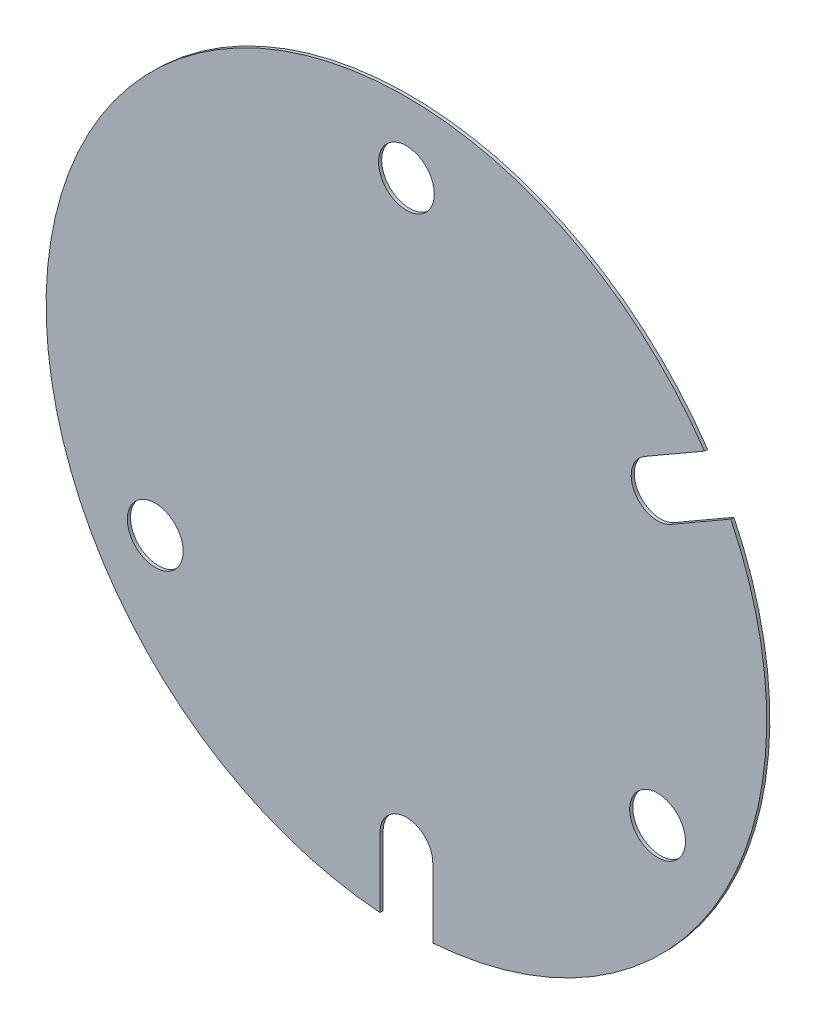
SolidWorks part; units mm, degrees
material "Copper"
ref_plane "Front Plane" through (0, 0, 0) normal (0, 0, 1) x (1, 0, 0)
ref_plane "Top Plane" through (0, 0, 0) normal (0, 1, 0) x (1, 0, 0)
ref_plane "Right Plane" through (0, 0, 0) normal (1, 0, 0) x (0, 0, -1)
sketch "Sketch3" plane through (0, 0, 0) normal (0, 0, 1) x (1, 0, 0)
  line L0 (0, 0) -> (0, 16.5) construction
  circle A0 centre (0, 0) radius 20.5
  circle A1 centre (0, 16.5) radius 1.5875
  circle A2 centre (14.2894, -8.25) radius 1.5875
  circle A3 centre (-14.2894, -8.25) radius 1.5875
  circle A4 centre (0, 0) radius 16.5 construction
  circle A6 centre (14.2894, -8.25) radius 1.5875
  circle A8 centre (-14.2894, -8.25) radius 1.5875
  circle A10 centre (-14.2894, 8.25) radius 1.5875 [skipped]
  circle A11 centre (0, -16.5) radius 1.5875 [skipped]
  circle A12 centre (14.2894, 8.25) radius 1.5875 [skipped]
  dimension "D1" = 41
  dimension "D2" = 3.175
  dimension "D3" = 33
  dimension "D4" = 3
  dimension "D5" = 6
extrude "Extrude2" add sketch "Sketch3" along normal blind 0.1778
sketch "Sketch5" plane through (0, 0, 0) normal (0, 0, 1) x (1, 0, 0)
  line L0 (1.5, -16.5) -> (1.5, -20.445)
  line L1 (-1.5, -16.5) -> (-1.5, -20.445)
  circle A0 centre (0, 0) radius 16.5 construction
  circle A1 centre (0, -16.5) radius 1.5
  dimension "D1" = 3
extrude "Cut-Extrude1" cut sketch "Sketch5" along normal through all
ref_axis "Axis1" through (0, 0, 0.1778) along (0, 0, -1)
pattern_circular "CirPattern1" count 3 over 360 about axis through (0, 0, 0.1778) along (0, 0, -1) skipping 1 of "Cut-Extrude1"
sketch "Sketch7" plane through (0, 0, 0.1778) normal (0, 0, 1) x (1, 0, 0)
  line L6 (18.4559, 8.9235) -> (15.0394, 6.951)
  line L7 (13.5394, 9.549) -> (16.9559, 11.5216)
  line L10 (-1.5, -20.445) -> (-1.5, -16.5)
  line L11 (1.5, -16.5) -> (1.5, -20.445)
  line L12 (18.4559, 8.9235) -> (15.0394, 6.951)
  line L13 (13.5394, 9.549) -> (16.9559, 11.5216)
  line L16 (-1.5, -20.445) -> (-1.5, -16.5)
  line L17 (1.5, -16.5) -> (1.5, -20.445)
  circle A0 centre (-14.2894, -8.25) radius 1.5875 construction
  circle A1 centre (0, 16.5) radius 1.5875 construction
  circle A2 centre (14.2894, -8.25) radius 1.5875 construction
  circle A3 centre (-14.2894, -8.25) radius 1.5875
  circle A4 centre (0, 16.5) radius 1.5875
  circle A5 centre (14.2894, -8.25) radius 1.5875
  arc A6 (1.5, -20.445) -> (18.4559, 8.9235) centre (0, 0) ccw
  arc A7 (13.5394, 9.549) -> (15.0394, 6.951) centre (14.2894, 8.25) ccw
  arc A8 (16.9559, 11.5216) -> (-1.5, -20.445) centre (0, 0) ccw
  arc A11 (1.5, -16.5) -> (-1.5, -16.5) centre (0, -16.5) ccw
  arc A12 (1.5, -20.445) -> (18.4559, 8.9235) centre (0, 0) ccw
  arc A13 (13.5394, 9.549) -> (15.0394, 6.951) centre (14.2894, 8.25) ccw
  arc A14 (16.9559, 11.5216) -> (-1.5, -20.445) centre (0, 0) ccw
  arc A17 (1.5, -16.5) -> (-1.5, -16.5) centre (0, -16.5) ccw
  dimension "D1" = 0
sketch "Sketch6" plane through (0, 0, 0.1778) normal (0, 0, 1) x (1, 0, 0)
  line L0 (0, 13.5) -> (0, 0)
  line L1 (0.5, 0) -> (0.25, 0.433)
  line L2 (0.25, 0.433) -> (-0.25, 0.433)
  line L3 (-0.25, 0.433) -> (-0.5, 0)
  line L4 (-0.5, 0) -> (-0.25, -0.433)
  line L5 (-0.25, -0.433) -> (0.25, -0.433)
  line L6 (0.25, -0.433) -> (0.5, 0)
  line L7 (1.382, 0.5092) -> (1.132, 0.9422)
  line L8 (1.132, 0.9422) -> (0.632, 0.9422)
  line L9 (0.632, 0.9422) -> (0.382, 0.5092)
  line L10 (0.382, 0.5092) -> (0.632, 0.0762)
  line L11 (0.632, 0.0762) -> (1.132, 0.0762)
  line L12 (1.132, 0.0762) -> (1.382, 0.5092)
  line L13 (0, 0) -> (13.5, 0)
  line L14 (2.01, 0.433) -> (1.51, 0.433)
  line L15 (1.51, 0.433) -> (1.26, 0)
  line L16 (1.26, 0) -> (1.51, -0.433)
  line L17 (1.51, -0.433) -> (2.01, -0.433)
  line L18 (2.01, -0.433) -> (2.26, 0)
  line L19 (2.26, 0) -> (2.01, 0.433)
  line L20 (2.142, 0.5092) -> (2.392, 0.0762)
  line L21 (2.392, 0.9422) -> (2.142, 0.5092)
  line L22 (2.892, 0.9422) -> (2.392, 0.9422)
  line L23 (3.142, 0.5092) -> (2.892, 0.9422)
  line L24 (2.892, 0.0762) -> (3.142, 0.5092)
  line L25 (2.392, 0.0762) -> (2.892, 0.0762)
  line L26 (3.77, 0.433) -> (3.27, 0.433)
  line L27 (3.27, 0.433) -> (3.02, 0)
  line L28 (3.02, 0) -> (3.27, -0.433)
  line L29 (3.27, -0.433) -> (3.77, -0.433)
  line L30 (3.77, -0.433) -> (4.02, 0)
  line L31 (4.02, 0) -> (3.77, 0.433)
  line L32 (3.902, 0.5092) -> (4.152, 0.0762)
  line L33 (4.152, 0.9422) -> (3.902, 0.5092)
  line L34 (4.652, 0.9422) -> (4.152, 0.9422)
  line L35 (4.902, 0.5092) -> (4.652, 0.9422)
  line L36 (4.652, 0.0762) -> (4.902, 0.5092)
  line L37 (4.152, 0.0762) -> (4.652, 0.0762)
  line L38 (5.53, 0.433) -> (5.03, 0.433)
  line L39 (5.03, 0.433) -> (4.78, 0)
  line L40 (4.78, 0) -> (5.03, -0.433)
  line L41 (5.03, -0.433) -> (5.53, -0.433)
  line L42 (5.53, -0.433) -> (5.78, 0)
  line L43 (5.78, 0) -> (5.53, 0.433)
  line L44 (5.662, 0.5092) -> (5.912, 0.0762)
  line L45 (5.912, 0.9422) -> (5.662, 0.5092)
  line L46 (6.412, 0.9422) -> (5.912, 0.9422)
  line L47 (6.662, 0.5092) -> (6.412, 0.9422)
  line L48 (6.412, 0.0762) -> (6.662, 0.5092)
  line L49 (5.912, 0.0762) -> (6.412, 0.0762)
  line L50 (7.29, 0.433) -> (6.79, 0.433)
  line L51 (6.79, 0.433) -> (6.54, 0)
  line L52 (6.54, 0) -> (6.79, -0.433)
  line L53 (6.79, -0.433) -> (7.29, -0.433)
  line L54 (7.29, -0.433) -> (7.54, 0)
  line L55 (7.54, 0) -> (7.29, 0.433)
  line L56 (7.422, 0.5092) -> (7.672, 0.0762)
  line L57 (7.672, 0.9422) -> (7.422, 0.5092)
  line L58 (8.172, 0.9422) -> (7.672, 0.9422)
  line L59 (8.422, 0.5092) -> (8.172, 0.9422)
  line L60 (8.172, 0.0762) -> (8.422, 0.5092)
  line L61 (7.672, 0.0762) -> (8.172, 0.0762)
  line L62 (9.05, 0.433) -> (8.55, 0.433)
  line L63 (8.55, 0.433) -> (8.3, 0)
  line L64 (8.3, 0) -> (8.55, -0.433)
  line L65 (8.55, -0.433) -> (9.05, -0.433)
  line L66 (9.05, -0.433) -> (9.3, 0)
  line L67 (9.3, 0) -> (9.05, 0.433)
  line L68 (9.182, 0.5092) -> (9.432, 0.0762)
  line L69 (9.432, 0.9422) -> (9.182, 0.5092)
  line L70 (9.932, 0.9422) -> (9.432, 0.9422)
  line L71 (10.182, 0.5092) -> (9.932, 0.9422)
  line L72 (9.932, 0.0762) -> (10.182, 0.5092)
  line L73 (9.432, 0.0762) -> (9.932, 0.0762)
  line L74 (10.81, 0.433) -> (10.31, 0.433)
  line L75 (10.31, 0.433) -> (10.06, 0)
  line L76 (10.06, 0) -> (10.31, -0.433)
  line L77 (10.31, -0.433) -> (10.81, -0.433)
  line L78 (10.81, -0.433) -> (11.06, 0)
  line L79 (11.06, 0) -> (10.81, 0.433)
  line L80 (10.942, 0.5092) -> (11.192, 0.0762)
  line L81 (11.192, 0.9422) -> (10.942, 0.5092)
  line L82 (11.692, 0.9422) -> (11.192, 0.9422)
  line L83 (11.942, 0.5092) -> (11.692, 0.9422)
  line L84 (11.692, 0.0762) -> (11.942, 0.5092)
  line L85 (11.192, 0.0762) -> (11.692, 0.0762)
  line L86 (12.57, 0.433) -> (12.07, 0.433)
  line L87 (12.07, 0.433) -> (11.82, 0)
  line L88 (11.82, 0) -> (12.07, -0.433)
  line L89 (12.07, -0.433) -> (12.57, -0.433)
  line L90 (12.57, -0.433) -> (12.82, 0)
  line L91 (12.82, 0) -> (12.57, 0.433)
  line L92 (12.702, 0.5092) -> (12.952, 0.0762)
  line L93 (12.952, 0.9422) -> (12.702, 0.5092)
  line L94 (13.452, 0.9422) -> (12.952, 0.9422)
  line L95 (13.702, 0.5092) -> (13.452, 0.9422)
  line L96 (13.452, 0.0762) -> (13.702, 0.5092)
  line L97 (12.952, 0.0762) -> (13.452, 0.0762)
  line L98 (14.33, 0.433) -> (13.83, 0.433)
  line L99 (13.83, 0.433) -> (13.58, 0)
  line L100 (13.58, 0) -> (13.83, -0.433)
  line L101 (13.83, -0.433) -> (14.33, -0.433)
  line L102 (14.33, -0.433) -> (14.58, 0)
  line L103 (14.58, 0) -> (14.33, 0.433)
  line L104 (14.462, 0.5092) -> (14.712, 0.0762)
  line L105 (14.712, 0.9422) -> (14.462, 0.5092)
  line L106 (15.212, 0.9422) -> (14.712, 0.9422)
  line L107 (15.462, 0.5092) -> (15.212, 0.9422)
  line L108 (15.212, 0.0762) -> (15.462, 0.5092)
  line L109 (14.712, 0.0762) -> (15.212, 0.0762)
  line L110 (0.25, 1.453) -> (-0.25, 1.453)
  line L111 (-0.25, 1.453) -> (-0.5, 1.02)
  line L112 (-0.5, 1.02) -> (-0.25, 0.587)
  line L113 (-0.25, 0.587) -> (0.25, 0.587)
  line L114 (0.25, 0.587) -> (0.5, 1.02)
  line L115 (0.5, 1.02) -> (0.25, 1.453)
  line L116 (0.382, 1.5292) -> (0.632, 1.0962)
  line L117 (0.632, 1.9622) -> (0.382, 1.5292)
  line L118 (1.132, 1.9622) -> (0.632, 1.9622)
  line L119 (1.382, 1.5292) -> (1.132, 1.9622)
  line L120 (1.132, 1.0962) -> (1.382, 1.5292)
  line L121 (0.632, 1.0962) -> (1.132, 1.0962)
  line L122 (2.01, 1.453) -> (1.51, 1.453)
  line L123 (1.51, 1.453) -> (1.26, 1.02)
  line L124 (1.26, 1.02) -> (1.51, 0.587)
  line L125 (1.51, 0.587) -> (2.01, 0.587)
  line L126 (2.01, 0.587) -> (2.26, 1.02)
  line L127 (2.26, 1.02) -> (2.01, 1.453)
  line L128 (2.142, 1.5292) -> (2.392, 1.0962)
  line L129 (2.392, 1.9622) -> (2.142, 1.5292)
  line L130 (2.892, 1.9622) -> (2.392, 1.9622)
  line L131 (3.142, 1.5292) -> (2.892, 1.9622)
  line L132 (2.892, 1.0962) -> (3.142, 1.5292)
  line L133 (2.392, 1.0962) -> (2.892, 1.0962)
  line L134 (3.77, 1.453) -> (3.27, 1.453)
  line L135 (3.27, 1.453) -> (3.02, 1.02)
  line L136 (3.02, 1.02) -> (3.27, 0.587)
  line L137 (3.27, 0.587) -> (3.77, 0.587)
  line L138 (3.77, 0.587) -> (4.02, 1.02)
  line L139 (4.02, 1.02) -> (3.77, 1.453)
  line L140 (3.902, 1.5292) -> (4.152, 1.0962)
  line L141 (4.152, 1.9622) -> (3.902, 1.5292)
  line L142 (4.652, 1.9622) -> (4.152, 1.9622)
  line L143 (4.902, 1.5292) -> (4.652, 1.9622)
  line L144 (4.652, 1.0962) -> (4.902, 1.5292)
  line L145 (4.152, 1.0962) -> (4.652, 1.0962)
  line L146 (5.53, 1.453) -> (5.03, 1.453)
  line L147 (5.03, 1.453) -> (4.78, 1.02)
  line L148 (4.78, 1.02) -> (5.03, 0.587)
  line L149 (5.03, 0.587) -> (5.53, 0.587)
  line L150 (5.53, 0.587) -> (5.78, 1.02)
  line L151 (5.78, 1.02) -> (5.53, 1.453)
  line L152 (5.662, 1.5292) -> (5.912, 1.0962)
  line L153 (5.912, 1.9622) -> (5.662, 1.5292)
  line L154 (6.412, 1.9622) -> (5.912, 1.9622)
  line L155 (6.662, 1.5292) -> (6.412, 1.9622)
  line L156 (6.412, 1.0962) -> (6.662, 1.5292)
  line L157 (5.912, 1.0962) -> (6.412, 1.0962)
  line L158 (7.29, 1.453) -> (6.79, 1.453)
  line L159 (6.79, 1.453) -> (6.54, 1.02)
  line L160 (6.54, 1.02) -> (6.79, 0.587)
  line L161 (6.79, 0.587) -> (7.29, 0.587)
  line L162 (7.29, 0.587) -> (7.54, 1.02)
  line L163 (7.54, 1.02) -> (7.29, 1.453)
  line L164 (7.422, 1.5292) -> (7.672, 1.0962)
  line L165 (7.672, 1.9622) -> (7.422, 1.5292)
  line L166 (8.172, 1.9622) -> (7.672, 1.9622)
  line L167 (8.422, 1.5292) -> (8.172, 1.9622)
  line L168 (8.172, 1.0962) -> (8.422, 1.5292)
  line L169 (7.672, 1.0962) -> (8.172, 1.0962)
  line L170 (9.05, 1.453) -> (8.55, 1.453)
  line L171 (8.55, 1.453) -> (8.3, 1.02)
  line L172 (8.3, 1.02) -> (8.55, 0.587)
  line L173 (8.55, 0.587) -> (9.05, 0.587)
  line L174 (9.05, 0.587) -> (9.3, 1.02)
  line L175 (9.3, 1.02) -> (9.05, 1.453)
  line L176 (9.182, 1.5292) -> (9.432, 1.0962)
  line L177 (9.432, 1.9622) -> (9.182, 1.5292)
  line L178 (9.932, 1.9622) -> (9.432, 1.9622)
  line L179 (10.182, 1.5292) -> (9.932, 1.9622)
  line L180 (9.932, 1.0962) -> (10.182, 1.5292)
  line L181 (9.432, 1.0962) -> (9.932, 1.0962)
  line L182 (10.81, 1.453) -> (10.31, 1.453)
  line L183 (10.31, 1.453) -> (10.06, 1.02)
  line L184 (10.06, 1.02) -> (10.31, 0.587)
  line L185 (10.31, 0.587) -> (10.81, 0.587)
  line L186 (10.81, 0.587) -> (11.06, 1.02)
  line L187 (11.06, 1.02) -> (10.81, 1.453)
  line L188 (10.942, 1.5292) -> (11.192, 1.0962)
  line L189 (11.192, 1.9622) -> (10.942, 1.5292)
  line L190 (11.692, 1.9622) -> (11.192, 1.9622)
  line L191 (11.942, 1.5292) -> (11.692, 1.9622)
  line L192 (11.692, 1.0962) -> (11.942, 1.5292)
  line L193 (11.192, 1.0962) -> (11.692, 1.0962)
  line L194 (12.57, 1.453) -> (12.07, 1.453)
  line L195 (12.07, 1.453) -> (11.82, 1.02)
  line L196 (11.82, 1.02) -> (12.07, 0.587)
  line L197 (12.07, 0.587) -> (12.57, 0.587)
  line L198 (12.57, 0.587) -> (12.82, 1.02)
  line L199 (12.82, 1.02) -> (12.57, 1.453)
  line L200 (12.702, 1.5292) -> (12.952, 1.0962)
  line L201 (12.952, 1.9622) -> (12.702, 1.5292)
  line L202 (13.452, 1.9622) -> (12.952, 1.9622)
  line L203 (13.702, 1.5292) -> (13.452, 1.9622)
  line L204 (13.452, 1.0962) -> (13.702, 1.5292)
  line L205 (12.952, 1.0962) -> (13.452, 1.0962)
  line L206 (14.33, 1.453) -> (13.83, 1.453)
  line L207 (13.83, 1.453) -> (13.58, 1.02)
  line L208 (13.58, 1.02) -> (13.83, 0.587)
  line L209 (13.83, 0.587) -> (14.33, 0.587)
  line L210 (14.33, 0.587) -> (14.58, 1.02)
  line L211 (14.58, 1.02) -> (14.33, 1.453)
  line L212 (14.462, 1.5292) -> (14.712, 1.0962)
  line L213 (14.712, 1.9622) -> (14.462, 1.5292)
  line L214 (15.212, 1.9622) -> (14.712, 1.9622)
  line L215 (15.462, 1.5292) -> (15.212, 1.9622)
  line L216 (15.212, 1.0962) -> (15.462, 1.5292)
  line L217 (14.712, 1.0962) -> (15.212, 1.0962)
  line L218 (0.25, 2.473) -> (-0.25, 2.473)
  line L219 (-0.25, 2.473) -> (-0.5, 2.04)
  line L220 (-0.5, 2.04) -> (-0.25, 1.607)
  line L221 (-0.25, 1.607) -> (0.25, 1.607)
  line L222 (0.25, 1.607) -> (0.5, 2.04)
  line L223 (0.5, 2.04) -> (0.25, 2.473)
  line L224 (0.382, 2.5492) -> (0.632, 2.1162)
  line L225 (0.632, 2.9822) -> (0.382, 2.5492)
  line L226 (1.132, 2.9822) -> (0.632, 2.9822)
  line L227 (1.382, 2.5492) -> (1.132, 2.9822)
  line L228 (1.132, 2.1162) -> (1.382, 2.5492)
  line L229 (0.632, 2.1162) -> (1.132, 2.1162)
  line L230 (2.01, 2.473) -> (1.51, 2.473)
  line L231 (1.51, 2.473) -> (1.26, 2.04)
  line L232 (1.26, 2.04) -> (1.51, 1.607)
  line L233 (1.51, 1.607) -> (2.01, 1.607)
  line L234 (2.01, 1.607) -> (2.26, 2.04)
  line L235 (2.26, 2.04) -> (2.01, 2.473)
  line L236 (2.142, 2.5492) -> (2.392, 2.1162)
  line L237 (2.392, 2.9822) -> (2.142, 2.5492)
  line L238 (2.892, 2.9822) -> (2.392, 2.9822)
  line L239 (3.142, 2.5492) -> (2.892, 2.9822)
  line L240 (2.892, 2.1162) -> (3.142, 2.5492)
  line L241 (2.392, 2.1162) -> (2.892, 2.1162)
  line L242 (3.77, 2.473) -> (3.27, 2.473)
  line L243 (3.27, 2.473) -> (3.02, 2.04)
  line L244 (3.02, 2.04) -> (3.27, 1.607)
  line L245 (3.27, 1.607) -> (3.77, 1.607)
  line L246 (3.77, 1.607) -> (4.02, 2.04)
  line L247 (4.02, 2.04) -> (3.77, 2.473)
  line L248 (3.902, 2.5492) -> (4.152, 2.1162)
  line L249 (4.152, 2.9822) -> (3.902, 2.5492)
  line L250 (4.652, 2.9822) -> (4.152, 2.9822)
  line L251 (4.902, 2.5492) -> (4.652, 2.9822)
  line L252 (4.652, 2.1162) -> (4.902, 2.5492)
  line L253 (4.152, 2.1162) -> (4.652, 2.1162)
  line L254 (5.53, 2.473) -> (5.03, 2.473)
  line L255 (5.03, 2.473) -> (4.78, 2.04)
  line L256 (4.78, 2.04) -> (5.03, 1.607)
  line L257 (5.03, 1.607) -> (5.53, 1.607)
  line L258 (5.53, 1.607) -> (5.78, 2.04)
  line L259 (5.78, 2.04) -> (5.53, 2.473)
  line L260 (5.662, 2.5492) -> (5.912, 2.1162)
  line L261 (5.912, 2.9822) -> (5.662, 2.5492)
  line L262 (6.412, 2.9822) -> (5.912, 2.9822)
  line L263 (6.662, 2.5492) -> (6.412, 2.9822)
  line L264 (6.412, 2.1162) -> (6.662, 2.5492)
  line L265 (5.912, 2.1162) -> (6.412, 2.1162)
  line L266 (7.29, 2.473) -> (6.79, 2.473)
  line L267 (6.79, 2.473) -> (6.54, 2.04)
  line L268 (6.54, 2.04) -> (6.79, 1.607)
  line L269 (6.79, 1.607) -> (7.29, 1.607)
  line L270 (7.29, 1.607) -> (7.54, 2.04)
  line L271 (7.54, 2.04) -> (7.29, 2.473)
  line L272 (7.422, 2.5492) -> (7.672, 2.1162)
  line L273 (7.672, 2.9822) -> (7.422, 2.5492)
  line L274 (8.172, 2.9822) -> (7.672, 2.9822)
  line L275 (8.422, 2.5492) -> (8.172, 2.9822)
  line L276 (8.172, 2.1162) -> (8.422, 2.5492)
  line L277 (7.672, 2.1162) -> (8.172, 2.1162)
  line L278 (9.05, 2.473) -> (8.55, 2.473)
  line L279 (8.55, 2.473) -> (8.3, 2.04)
  line L280 (8.3, 2.04) -> (8.55, 1.607)
  line L281 (8.55, 1.607) -> (9.05, 1.607)
  line L282 (9.05, 1.607) -> (9.3, 2.04)
  line L283 (9.3, 2.04) -> (9.05, 2.473)
  line L284 (9.182, 2.5492) -> (9.432, 2.1162)
  line L285 (9.432, 2.9822) -> (9.182, 2.5492)
  line L286 (9.932, 2.9822) -> (9.432, 2.9822)
  line L287 (10.182, 2.5492) -> (9.932, 2.9822)
  line L288 (9.932, 2.1162) -> (10.182, 2.5492)
  line L289 (9.432, 2.1162) -> (9.932, 2.1162)
  line L290 (10.81, 2.473) -> (10.31, 2.473)
  line L291 (10.31, 2.473) -> (10.06, 2.04)
  line L292 (10.06, 2.04) -> (10.31, 1.607)
  line L293 (10.31, 1.607) -> (10.81, 1.607)
  line L294 (10.81, 1.607) -> (11.06, 2.04)
  line L295 (11.06, 2.04) -> (10.81, 2.473)
  line L296 (10.942, 2.5492) -> (11.192, 2.1162)
  line L297 (11.192, 2.9822) -> (10.942, 2.5492)
  line L298 (11.692, 2.9822) -> (11.192, 2.9822)
  line L299 (11.942, 2.5492) -> (11.692, 2.9822)
  line L300 (11.692, 2.1162) -> (11.942, 2.5492)
  line L301 (11.192, 2.1162) -> (11.692, 2.1162)
  line L302 (12.57, 2.473) -> (12.07, 2.473)
  line L303 (12.07, 2.473) -> (11.82, 2.04)
  line L304 (11.82, 2.04) -> (12.07, 1.607)
  line L305 (12.07, 1.607) -> (12.57, 1.607)
  line L306 (12.57, 1.607) -> (12.82, 2.04)
  line L307 (12.82, 2.04) -> (12.57, 2.473)
  line L308 (12.702, 2.5492) -> (12.952, 2.1162)
  line L309 (12.952, 2.9822) -> (12.702, 2.5492)
  line L310 (13.452, 2.9822) -> (12.952, 2.9822)
  line L311 (13.702, 2.5492) -> (13.452, 2.9822)
  line L312 (13.452, 2.1162) -> (13.702, 2.5492)
  line L313 (12.952, 2.1162) -> (13.452, 2.1162)
  line L314 (14.33, 2.473) -> (13.83, 2.473)
  line L315 (13.83, 2.473) -> (13.58, 2.04)
  line L316 (13.58, 2.04) -> (13.83, 1.607)
  line L317 (13.83, 1.607) -> (14.33, 1.607)
  line L318 (14.33, 1.607) -> (14.58, 2.04)
  line L319 (14.58, 2.04) -> (14.33, 2.473)
  line L320 (14.462, 2.5492) -> (14.712, 2.1162)
  line L321 (14.712, 2.9822) -> (14.462, 2.5492)
  line L322 (15.212, 2.9822) -> (14.712, 2.9822)
  line L323 (15.462, 2.5492) -> (15.212, 2.9822)
  line L324 (15.212, 2.1162) -> (15.462, 2.5492)
  line L325 (14.712, 2.1162) -> (15.212, 2.1162)
  line L326 (0.25, 3.493) -> (-0.25, 3.493)
  line L327 (-0.25, 3.493) -> (-0.5, 3.06)
  line L328 (-0.5, 3.06) -> (-0.25, 2.627)
  line L329 (-0.25, 2.627) -> (0.25, 2.627)
  line L330 (0.25, 2.627) -> (0.5, 3.06)
  line L331 (0.5, 3.06) -> (0.25, 3.493)
  line L332 (0.382, 3.5692) -> (0.632, 3.1362)
  line L333 (0.632, 4.0022) -> (0.382, 3.5692)
  line L334 (1.132, 4.0022) -> (0.632, 4.0022)
  line L335 (1.382, 3.5692) -> (1.132, 4.0022)
  line L336 (1.132, 3.1362) -> (1.382, 3.5692)
  line L337 (0.632, 3.1362) -> (1.132, 3.1362)
  line L338 (2.01, 3.493) -> (1.51, 3.493)
  line L339 (1.51, 3.493) -> (1.26, 3.06)
  line L340 (1.26, 3.06) -> (1.51, 2.627)
  line L341 (1.51, 2.627) -> (2.01, 2.627)
  line L342 (2.01, 2.627) -> (2.26, 3.06)
  line L343 (2.26, 3.06) -> (2.01, 3.493)
  line L344 (2.142, 3.5692) -> (2.392, 3.1362)
  line L345 (2.392, 4.0022) -> (2.142, 3.5692)
  line L346 (2.892, 4.0022) -> (2.392, 4.0022)
  line L347 (3.142, 3.5692) -> (2.892, 4.0022)
  line L348 (2.892, 3.1362) -> (3.142, 3.5692)
  line L349 (2.392, 3.1362) -> (2.892, 3.1362)
  line L350 (3.77, 3.493) -> (3.27, 3.493)
  line L351 (3.27, 3.493) -> (3.02, 3.06)
  line L352 (3.02, 3.06) -> (3.27, 2.627)
  line L353 (3.27, 2.627) -> (3.77, 2.627)
  line L354 (3.77, 2.627) -> (4.02, 3.06)
  line L355 (4.02, 3.06) -> (3.77, 3.493)
  line L356 (3.902, 3.5692) -> (4.152, 3.1362)
  line L357 (4.152, 4.0022) -> (3.902, 3.5692)
  line L358 (4.652, 4.0022) -> (4.152, 4.0022)
  line L359 (4.902, 3.5692) -> (4.652, 4.0022)
  line L360 (4.652, 3.1362) -> (4.902, 3.5692)
  line L361 (4.152, 3.1362) -> (4.652, 3.1362)
  line L362 (5.53, 3.493) -> (5.03, 3.493)
  line L363 (5.03, 3.493) -> (4.78, 3.06)
  line L364 (4.78, 3.06) -> (5.03, 2.627)
  line L365 (5.03, 2.627) -> (5.53, 2.627)
  line L366 (5.53, 2.627) -> (5.78, 3.06)
  line L367 (5.78, 3.06) -> (5.53, 3.493)
  line L368 (5.662, 3.5692) -> (5.912, 3.1362)
  line L369 (5.912, 4.0022) -> (5.662, 3.5692)
  line L370 (6.412, 4.0022) -> (5.912, 4.0022)
  line L371 (6.662, 3.5692) -> (6.412, 4.0022)
  line L372 (6.412, 3.1362) -> (6.662, 3.5692)
  line L373 (5.912, 3.1362) -> (6.412, 3.1362)
  line L374 (7.29, 3.493) -> (6.79, 3.493)
  line L375 (6.79, 3.493) -> (6.54, 3.06)
  line L376 (6.54, 3.06) -> (6.79, 2.627)
  line L377 (6.79, 2.627) -> (7.29, 2.627)
  line L378 (7.29, 2.627) -> (7.54, 3.06)
  line L379 (7.54, 3.06) -> (7.29, 3.493)
  line L380 (7.422, 3.5692) -> (7.672, 3.1362)
  line L381 (7.672, 4.0022) -> (7.422, 3.5692)
  line L382 (8.172, 4.0022) -> (7.672, 4.0022)
  line L383 (8.422, 3.5692) -> (8.172, 4.0022)
  line L384 (8.172, 3.1362) -> (8.422, 3.5692)
  line L385 (7.672, 3.1362) -> (8.172, 3.1362)
  line L386 (9.05, 3.493) -> (8.55, 3.493)
  line L387 (8.55, 3.493) -> (8.3, 3.06)
  line L388 (8.3, 3.06) -> (8.55, 2.627)
  line L389 (8.55, 2.627) -> (9.05, 2.627)
  line L390 (9.05, 2.627) -> (9.3, 3.06)
  line L391 (9.3, 3.06) -> (9.05, 3.493)
  line L392 (9.182, 3.5692) -> (9.432, 3.1362)
  line L393 (9.432, 4.0022) -> (9.182, 3.5692)
  line L394 (9.932, 4.0022) -> (9.432, 4.0022)
  line L395 (10.182, 3.5692) -> (9.932, 4.0022)
  line L396 (9.932, 3.1362) -> (10.182, 3.5692)
  line L397 (9.432, 3.1362) -> (9.932, 3.1362)
  line L398 (10.81, 3.493) -> (10.31, 3.493)
  line L399 (10.31, 3.493) -> (10.06, 3.06)
  line L400 (10.06, 3.06) -> (10.31, 2.627)
  line L401 (10.31, 2.627) -> (10.81, 2.627)
  line L402 (10.81, 2.627) -> (11.06, 3.06)
  line L403 (11.06, 3.06) -> (10.81, 3.493)
  line L404 (10.942, 3.5692) -> (11.192, 3.1362)
  line L405 (11.192, 4.0022) -> (10.942, 3.5692)
  line L406 (11.692, 4.0022) -> (11.192, 4.0022)
  line L407 (11.942, 3.5692) -> (11.692, 4.0022)
  line L408 (11.692, 3.1362) -> (11.942, 3.5692)
  line L409 (11.192, 3.1362) -> (11.692, 3.1362)
  line L410 (12.57, 3.493) -> (12.07, 3.493)
  line L411 (12.07, 3.493) -> (11.82, 3.06)
  line L412 (11.82, 3.06) -> (12.07, 2.627)
  line L413 (12.07, 2.627) -> (12.57, 2.627)
  line L414 (12.57, 2.627) -> (12.82, 3.06)
  line L415 (12.82, 3.06) -> (12.57, 3.493)
  line L416 (12.702, 3.5692) -> (12.952, 3.1362)
  line L417 (12.952, 4.0022) -> (12.702, 3.5692)
  line L418 (13.452, 4.0022) -> (12.952, 4.0022)
  line L419 (13.702, 3.5692) -> (13.452, 4.0022)
  line L420 (13.452, 3.1362) -> (13.702, 3.5692)
  line L421 (12.952, 3.1362) -> (13.452, 3.1362)
  line L422 (14.33, 3.493) -> (13.83, 3.493)
  line L423 (13.83, 3.493) -> (13.58, 3.06)
  line L424 (13.58, 3.06) -> (13.83, 2.627)
  line L425 (13.83, 2.627) -> (14.33, 2.627)
  line L426 (14.33, 2.627) -> (14.58, 3.06)
  line L427 (14.58, 3.06) -> (14.33, 3.493)
  line L428 (14.462, 3.5692) -> (14.712, 3.1362)
  line L429 (14.712, 4.0022) -> (14.462, 3.5692)
  line L430 (15.212, 4.0022) -> (14.712, 4.0022)
  line L431 (15.462, 3.5692) -> (15.212, 4.0022)
  line L432 (15.212, 3.1362) -> (15.462, 3.5692)
  line L433 (14.712, 3.1362) -> (15.212, 3.1362)
  line L434 (0.25, 4.513) -> (-0.25, 4.513)
  line L435 (-0.25, 4.513) -> (-0.5, 4.08)
  line L436 (-0.5, 4.08) -> (-0.25, 3.647)
  line L437 (-0.25, 3.647) -> (0.25, 3.647)
  line L438 (0.25, 3.647) -> (0.5, 4.08)
  line L439 (0.5, 4.08) -> (0.25, 4.513)
  line L440 (0.382, 4.5892) -> (0.632, 4.1562)
  line L441 (0.632, 5.0222) -> (0.382, 4.5892)
  line L442 (1.132, 5.0222) -> (0.632, 5.0222)
  line L443 (1.382, 4.5892) -> (1.132, 5.0222)
  line L444 (1.132, 4.1562) -> (1.382, 4.5892)
  line L445 (0.632, 4.1562) -> (1.132, 4.1562)
  line L446 (2.01, 4.513) -> (1.51, 4.513)
  line L447 (1.51, 4.513) -> (1.26, 4.08)
  line L448 (1.26, 4.08) -> (1.51, 3.647)
  line L449 (1.51, 3.647) -> (2.01, 3.647)
  line L450 (2.01, 3.647) -> (2.26, 4.08)
  line L451 (2.26, 4.08) -> (2.01, 4.513)
  line L452 (2.142, 4.5892) -> (2.392, 4.1562)
  line L453 (2.392, 5.0222) -> (2.142, 4.5892)
  line L454 (2.892, 5.0222) -> (2.392, 5.0222)
  line L455 (3.142, 4.5892) -> (2.892, 5.0222)
  line L456 (2.892, 4.1562) -> (3.142, 4.5892)
  line L457 (2.392, 4.1562) -> (2.892, 4.1562)
  line L458 (3.77, 4.513) -> (3.27, 4.513)
  line L459 (3.27, 4.513) -> (3.02, 4.08)
  line L460 (3.02, 4.08) -> (3.27, 3.647)
  line L461 (3.27, 3.647) -> (3.77, 3.647)
  line L462 (3.77, 3.647) -> (4.02, 4.08)
  line L463 (4.02, 4.08) -> (3.77, 4.513)
  line L464 (3.902, 4.5892) -> (4.152, 4.1562)
  line L465 (4.152, 5.0222) -> (3.902, 4.5892)
  line L466 (4.652, 5.0222) -> (4.152, 5.0222)
  line L467 (4.902, 4.5892) -> (4.652, 5.0222)
  line L468 (4.652, 4.1562) -> (4.902, 4.5892)
  line L469 (4.152, 4.1562) -> (4.652, 4.1562)
  line L470 (5.53, 4.513) -> (5.03, 4.513)
  line L471 (5.03, 4.513) -> (4.78, 4.08)
  line L472 (4.78, 4.08) -> (5.03, 3.647)
  line L473 (5.03, 3.647) -> (5.53, 3.647)
  line L474 (5.53, 3.647) -> (5.78, 4.08)
  line L475 (5.78, 4.08) -> (5.53, 4.513)
  line L476 (5.662, 4.5892) -> (5.912, 4.1562)
  line L477 (5.912, 5.0222) -> (5.662, 4.5892)
  line L478 (6.412, 5.0222) -> (5.912, 5.0222)
  line L479 (6.662, 4.5892) -> (6.412, 5.0222)
  line L480 (6.412, 4.1562) -> (6.662, 4.5892)
  line L481 (5.912, 4.1562) -> (6.412, 4.1562)
  line L482 (7.29, 4.513) -> (6.79, 4.513)
  line L483 (6.79, 4.513) -> (6.54, 4.08)
  line L484 (6.54, 4.08) -> (6.79, 3.647)
  line L485 (6.79, 3.647) -> (7.29, 3.647)
  line L486 (7.29, 3.647) -> (7.54, 4.08)
  line L487 (7.54, 4.08) -> (7.29, 4.513)
  line L488 (7.422, 4.5892) -> (7.672, 4.1562)
  line L489 (7.672, 5.0222) -> (7.422, 4.5892)
  line L490 (8.172, 5.0222) -> (7.672, 5.0222)
  line L491 (8.422, 4.5892) -> (8.172, 5.0222)
  line L492 (8.172, 4.1562) -> (8.422, 4.5892)
  line L493 (7.672, 4.1562) -> (8.172, 4.1562)
  line L494 (9.05, 4.513) -> (8.55, 4.513)
  line L495 (8.55, 4.513) -> (8.3, 4.08)
  line L496 (8.3, 4.08) -> (8.55, 3.647)
  line L497 (8.55, 3.647) -> (9.05, 3.647)
  line L498 (9.05, 3.647) -> (9.3, 4.08)
  line L499 (9.3, 4.08) -> (9.05, 4.513)
  line L500 (9.182, 4.5892) -> (9.432, 4.1562)
  line L501 (9.432, 5.0222) -> (9.182, 4.5892)
  line L502 (9.932, 5.0222) -> (9.432, 5.0222)
  line L503 (10.182, 4.5892) -> (9.932, 5.0222)
  line L504 (9.932, 4.1562) -> (10.182, 4.5892)
  line L505 (9.432, 4.1562) -> (9.932, 4.1562)
  line L506 (10.81, 4.513) -> (10.31, 4.513)
  line L507 (10.31, 4.513) -> (10.06, 4.08)
  line L508 (10.06, 4.08) -> (10.31, 3.647)
  line L509 (10.31, 3.647) -> (10.81, 3.647)
  line L510 (10.81, 3.647) -> (11.06, 4.08)
  line L511 (11.06, 4.08) -> (10.81, 4.513)
  line L512 (10.942, 4.5892) -> (11.192, 4.1562)
  line L513 (11.192, 5.0222) -> (10.942, 4.5892)
  line L514 (11.692, 5.0222) -> (11.192, 5.0222)
  line L515 (11.942, 4.5892) -> (11.692, 5.0222)
  line L516 (11.692, 4.1562) -> (11.942, 4.5892)
  line L517 (11.192, 4.1562) -> (11.692, 4.1562)
  line L518 (12.57, 4.513) -> (12.07, 4.513)
  line L519 (12.07, 4.513) -> (11.82, 4.08)
  line L520 (11.82, 4.08) -> (12.07, 3.647)
  line L521 (12.07, 3.647) -> (12.57, 3.647)
  line L522 (12.57, 3.647) -> (12.82, 4.08)
  line L523 (12.82, 4.08) -> (12.57, 4.513)
  line L524 (12.702, 4.5892) -> (12.952, 4.1562)
  line L525 (12.952, 5.0222) -> (12.702, 4.5892)
  line L526 (13.452, 5.0222) -> (12.952, 5.0222)
  line L527 (13.702, 4.5892) -> (13.452, 5.0222)
  line L528 (13.452, 4.1562) -> (13.702, 4.5892)
  line L529 (12.952, 4.1562) -> (13.452, 4.1562)
  line L530 (14.33, 4.513) -> (13.83, 4.513)
  line L531 (13.83, 4.513) -> (13.58, 4.08)
  line L532 (13.58, 4.08) -> (13.83, 3.647)
  line L533 (13.83, 3.647) -> (14.33, 3.647)
  line L534 (14.33, 3.647) -> (14.58, 4.08)
  line L535 (14.58, 4.08) -> (14.33, 4.513)
  line L536 (14.462, 4.5892) -> (14.712, 4.1562)
  line L537 (14.712, 5.0222) -> (14.462, 4.5892)
  line L538 (15.212, 5.0222) -> (14.712, 5.0222)
  line L539 (15.462, 4.5892) -> (15.212, 5.0222)
  line L540 (15.212, 4.1562) -> (15.462, 4.5892)
  line L541 (14.712, 4.1562) -> (15.212, 4.1562)
  line L542 (0.25, 5.533) -> (-0.25, 5.533)
  line L543 (-0.25, 5.533) -> (-0.5, 5.1)
  line L544 (-0.5, 5.1) -> (-0.25, 4.667)
  line L545 (-0.25, 4.667) -> (0.25, 4.667)
  line L546 (0.25, 4.667) -> (0.5, 5.1)
  line L547 (0.5, 5.1) -> (0.25, 5.533)
  line L548 (0.382, 5.6092) -> (0.632, 5.1762)
  line L549 (0.632, 6.0422) -> (0.382, 5.6092)
  line L550 (1.132, 6.0422) -> (0.632, 6.0422)
  line L551 (1.382, 5.6092) -> (1.132, 6.0422)
  line L552 (1.132, 5.1762) -> (1.382, 5.6092)
  line L553 (0.632, 5.1762) -> (1.132, 5.1762)
  line L554 (2.01, 5.533) -> (1.51, 5.533)
  line L555 (1.51, 5.533) -> (1.26, 5.1)
  line L556 (1.26, 5.1) -> (1.51, 4.667)
  line L557 (1.51, 4.667) -> (2.01, 4.667)
  line L558 (2.01, 4.667) -> (2.26, 5.1)
  line L559 (2.26, 5.1) -> (2.01, 5.533)
  line L560 (2.142, 5.6092) -> (2.392, 5.1762)
  line L561 (2.392, 6.0422) -> (2.142, 5.6092)
  line L562 (2.892, 6.0422) -> (2.392, 6.0422)
  line L563 (3.142, 5.6092) -> (2.892, 6.0422)
  line L564 (2.892, 5.1762) -> (3.142, 5.6092)
  line L565 (2.392, 5.1762) -> (2.892, 5.1762)
  line L566 (3.77, 5.533) -> (3.27, 5.533)
  line L567 (3.27, 5.533) -> (3.02, 5.1)
  line L568 (3.02, 5.1) -> (3.27, 4.667)
  line L569 (3.27, 4.667) -> (3.77, 4.667)
  line L570 (3.77, 4.667) -> (4.02, 5.1)
  line L571 (4.02, 5.1) -> (3.77, 5.533)
  line L572 (3.902, 5.6092) -> (4.152, 5.1762)
  line L573 (4.152, 6.0422) -> (3.902, 5.6092)
  line L574 (4.652, 6.0422) -> (4.152, 6.0422)
  line L575 (4.902, 5.6092) -> (4.652, 6.0422)
  line L576 (4.652, 5.1762) -> (4.902, 5.6092)
  line L577 (4.152, 5.1762) -> (4.652, 5.1762)
  line L578 (5.53, 5.533) -> (5.03, 5.533)
  line L579 (5.03, 5.533) -> (4.78, 5.1)
  line L580 (4.78, 5.1) -> (5.03, 4.667)
  line L581 (5.03, 4.667) -> (5.53, 4.667)
  line L582 (5.53, 4.667) -> (5.78, 5.1)
  line L583 (5.78, 5.1) -> (5.53, 5.533)
  line L584 (5.662, 5.6092) -> (5.912, 5.1762)
  line L585 (5.912, 6.0422) -> (5.662, 5.6092)
  line L586 (6.412, 6.0422) -> (5.912, 6.0422)
  line L587 (6.662, 5.6092) -> (6.412, 6.0422)
  line L588 (6.412, 5.1762) -> (6.662, 5.6092)
  line L589 (5.912, 5.1762) -> (6.412, 5.1762)
  line L590 (7.29, 5.533) -> (6.79, 5.533)
  line L591 (6.79, 5.533) -> (6.54, 5.1)
  line L592 (6.54, 5.1) -> (6.79, 4.667)
  line L593 (6.79, 4.667) -> (7.29, 4.667)
  line L594 (7.29, 4.667) -> (7.54, 5.1)
  line L595 (7.54, 5.1) -> (7.29, 5.533)
  line L596 (7.422, 5.6092) -> (7.672, 5.1762)
  line L597 (7.672, 6.0422) -> (7.422, 5.6092)
  line L598 (8.172, 6.0422) -> (7.672, 6.0422)
  line L599 (8.422, 5.6092) -> (8.172, 6.0422)
  line L600 (8.172, 5.1762) -> (8.422, 5.6092)
  line L601 (7.672, 5.1762) -> (8.172, 5.1762)
  line L602 (9.05, 5.533) -> (8.55, 5.533)
  line L603 (8.55, 5.533) -> (8.3, 5.1)
  line L604 (8.3, 5.1) -> (8.55, 4.667)
  line L605 (8.55, 4.667) -> (9.05, 4.667)
  line L606 (9.05, 4.667) -> (9.3, 5.1)
  line L607 (9.3, 5.1) -> (9.05, 5.533)
  line L608 (9.182, 5.6092) -> (9.432, 5.1762)
  line L609 (9.432, 6.0422) -> (9.182, 5.6092)
  line L610 (9.932, 6.0422) -> (9.432, 6.0422)
  line L611 (10.182, 5.6092) -> (9.932, 6.0422)
  line L612 (9.932, 5.1762) -> (10.182, 5.6092)
  line L613 (9.432, 5.1762) -> (9.932, 5.1762)
  line L614 (10.81, 5.533) -> (10.31, 5.533)
  line L615 (10.31, 5.533) -> (10.06, 5.1)
  line L616 (10.06, 5.1) -> (10.31, 4.667)
  line L617 (10.31, 4.667) -> (10.81, 4.667)
  line L618 (10.81, 4.667) -> (11.06, 5.1)
  line L619 (11.06, 5.1) -> (10.81, 5.533)
  line L620 (10.942, 5.6092) -> (11.192, 5.1762)
  line L621 (11.192, 6.0422) -> (10.942, 5.6092)
  line L622 (11.692, 6.0422) -> (11.192, 6.0422)
  line L623 (11.942, 5.6092) -> (11.692, 6.0422)
  line L624 (11.692, 5.1762) -> (11.942, 5.6092)
  line L625 (11.192, 5.1762) -> (11.692, 5.1762)
  line L626 (12.57, 5.533) -> (12.07, 5.533)
  line L627 (12.07, 5.533) -> (11.82, 5.1)
  line L628 (11.82, 5.1) -> (12.07, 4.667)
  line L629 (12.07, 4.667) -> (12.57, 4.667)
  line L630 (12.57, 4.667) -> (12.82, 5.1)
  line L631 (12.82, 5.1) -> (12.57, 5.533)
  line L632 (12.702, 5.6092) -> (12.952, 5.1762)
  line L633 (12.952, 6.0422) -> (12.702, 5.6092)
  line L634 (13.452, 6.0422) -> (12.952, 6.0422)
  line L635 (13.702, 5.6092) -> (13.452, 6.0422)
  line L636 (13.452, 5.1762) -> (13.702, 5.6092)
  line L637 (12.952, 5.1762) -> (13.452, 5.1762)
  line L638 (14.33, 5.533) -> (13.83, 5.533)
  line L639 (13.83, 5.533) -> (13.58, 5.1)
  line L640 (13.58, 5.1) -> (13.83, 4.667)
  line L641 (13.83, 4.667) -> (14.33, 4.667)
  line L642 (14.33, 4.667) -> (14.58, 5.1)
  line L643 (14.58, 5.1) -> (14.33, 5.533)
  line L644 (14.462, 5.6092) -> (14.712, 5.1762)
  line L645 (14.712, 6.0422) -> (14.462, 5.6092)
  line L646 (15.212, 6.0422) -> (14.712, 6.0422)
  line L647 (15.462, 5.6092) -> (15.212, 6.0422)
  line L648 (15.212, 5.1762) -> (15.462, 5.6092)
  line L649 (14.712, 5.1762) -> (15.212, 5.1762)
  line L650 (0.25, 6.553) -> (-0.25, 6.553)
  line L651 (-0.25, 6.553) -> (-0.5, 6.12)
  line L652 (-0.5, 6.12) -> (-0.25, 5.687)
  line L653 (-0.25, 5.687) -> (0.25, 5.687)
  line L654 (0.25, 5.687) -> (0.5, 6.12)
  line L655 (0.5, 6.12) -> (0.25, 6.553)
  line L656 (0.382, 6.6292) -> (0.632, 6.1962)
  line L657 (0.632, 7.0622) -> (0.382, 6.6292)
  line L658 (1.132, 7.0622) -> (0.632, 7.0622)
  line L659 (1.382, 6.6292) -> (1.132, 7.0622)
  line L660 (1.132, 6.1962) -> (1.382, 6.6292)
  line L661 (0.632, 6.1962) -> (1.132, 6.1962)
  line L662 (2.01, 6.553) -> (1.51, 6.553)
  line L663 (1.51, 6.553) -> (1.26, 6.12)
  line L664 (1.26, 6.12) -> (1.51, 5.687)
  line L665 (1.51, 5.687) -> (2.01, 5.687)
  line L666 (2.01, 5.687) -> (2.26, 6.12)
  line L667 (2.26, 6.12) -> (2.01, 6.553)
  line L668 (2.142, 6.6292) -> (2.392, 6.1962)
  line L669 (2.392, 7.0622) -> (2.142, 6.6292)
  line L670 (2.892, 7.0622) -> (2.392, 7.0622)
  line L671 (3.142, 6.6292) -> (2.892, 7.0622)
  line L672 (2.892, 6.1962) -> (3.142, 6.6292)
  line L673 (2.392, 6.1962) -> (2.892, 6.1962)
  line L674 (3.77, 6.553) -> (3.27, 6.553)
  line L675 (3.27, 6.553) -> (3.02, 6.12)
  line L676 (3.02, 6.12) -> (3.27, 5.687)
  line L677 (3.27, 5.687) -> (3.77, 5.687)
  line L678 (3.77, 5.687) -> (4.02, 6.12)
  line L679 (4.02, 6.12) -> (3.77, 6.553)
  line L680 (3.902, 6.6292) -> (4.152, 6.1962)
  line L681 (4.152, 7.0622) -> (3.902, 6.6292)
  line L682 (4.652, 7.0622) -> (4.152, 7.0622)
  line L683 (4.902, 6.6292) -> (4.652, 7.0622)
  line L684 (4.652, 6.1962) -> (4.902, 6.6292)
  line L685 (4.152, 6.1962) -> (4.652, 6.1962)
  line L686 (5.53, 6.553) -> (5.03, 6.553)
  line L687 (5.03, 6.553) -> (4.78, 6.12)
  line L688 (4.78, 6.12) -> (5.03, 5.687)
  line L689 (5.03, 5.687) -> (5.53, 5.687)
  line L690 (5.53, 5.687) -> (5.78, 6.12)
  line L691 (5.78, 6.12) -> (5.53, 6.553)
  line L692 (5.662, 6.6292) -> (5.912, 6.1962)
  line L693 (5.912, 7.0622) -> (5.662, 6.6292)
  line L694 (6.412, 7.0622) -> (5.912, 7.0622)
  line L695 (6.662, 6.6292) -> (6.412, 7.0622)
  line L696 (6.412, 6.1962) -> (6.662, 6.6292)
  line L697 (5.912, 6.1962) -> (6.412, 6.1962)
  line L698 (7.29, 6.553) -> (6.79, 6.553)
  line L699 (6.79, 6.553) -> (6.54, 6.12)
  line L700 (6.54, 6.12) -> (6.79, 5.687)
  line L701 (6.79, 5.687) -> (7.29, 5.687)
  line L702 (7.29, 5.687) -> (7.54, 6.12)
  line L703 (7.54, 6.12) -> (7.29, 6.553)
  line L704 (7.422, 6.6292) -> (7.672, 6.1962)
  line L705 (7.672, 7.0622) -> (7.422, 6.6292)
  line L706 (8.172, 7.0622) -> (7.672, 7.0622)
  line L707 (8.422, 6.6292) -> (8.172, 7.0622)
  line L708 (8.172, 6.1962) -> (8.422, 6.6292)
  line L709 (7.672, 6.1962) -> (8.172, 6.1962)
  line L710 (9.05, 6.553) -> (8.55, 6.553)
  line L711 (8.55, 6.553) -> (8.3, 6.12)
  line L712 (8.3, 6.12) -> (8.55, 5.687)
  line L713 (8.55, 5.687) -> (9.05, 5.687)
  line L714 (9.05, 5.687) -> (9.3, 6.12)
  line L715 (9.3, 6.12) -> (9.05, 6.553)
  line L716 (9.182, 6.6292) -> (9.432, 6.1962)
  line L717 (9.432, 7.0622) -> (9.182, 6.6292)
  line L718 (9.932, 7.0622) -> (9.432, 7.0622)
  line L719 (10.182, 6.6292) -> (9.932, 7.0622)
  line L720 (9.932, 6.1962) -> (10.182, 6.6292)
  line L721 (9.432, 6.1962) -> (9.932, 6.1962)
  line L722 (10.81, 6.553) -> (10.31, 6.553)
  line L723 (10.31, 6.553) -> (10.06, 6.12)
  line L724 (10.06, 6.12) -> (10.31, 5.687)
  line L725 (10.31, 5.687) -> (10.81, 5.687)
  line L726 (10.81, 5.687) -> (11.06, 6.12)
  line L727 (11.06, 6.12) -> (10.81, 6.553)
  line L728 (10.942, 6.6292) -> (11.192, 6.1962)
  line L729 (11.192, 7.0622) -> (10.942, 6.6292)
  line L730 (11.692, 7.0622) -> (11.192, 7.0622)
  line L731 (11.942, 6.6292) -> (11.692, 7.0622)
  line L732 (11.692, 6.1962) -> (11.942, 6.6292)
  line L733 (11.192, 6.1962) -> (11.692, 6.1962)
  line L734 (12.57, 6.553) -> (12.07, 6.553)
  line L735 (12.07, 6.553) -> (11.82, 6.12)
  line L736 (11.82, 6.12) -> (12.07, 5.687)
  line L737 (12.07, 5.687) -> (12.57, 5.687)
  line L738 (12.57, 5.687) -> (12.82, 6.12)
  line L739 (12.82, 6.12) -> (12.57, 6.553)
  line L740 (12.702, 6.6292) -> (12.952, 6.1962)
  line L741 (12.952, 7.0622) -> (12.702, 6.6292)
  line L742 (13.452, 7.0622) -> (12.952, 7.0622)
  line L743 (13.702, 6.6292) -> (13.452, 7.0622)
  line L744 (13.452, 6.1962) -> (13.702, 6.6292)
  line L745 (12.952, 6.1962) -> (13.452, 6.1962)
  line L746 (14.33, 6.553) -> (13.83, 6.553)
  line L747 (13.83, 6.553) -> (13.58, 6.12)
  line L748 (13.58, 6.12) -> (13.83, 5.687)
  line L749 (13.83, 5.687) -> (14.33, 5.687)
  line L750 (14.33, 5.687) -> (14.58, 6.12)
  line L751 (14.58, 6.12) -> (14.33, 6.553)
  line L752 (14.462, 6.6292) -> (14.712, 6.1962)
  line L753 (14.712, 7.0622) -> (14.462, 6.6292)
  line L754 (15.212, 7.0622) -> (14.712, 7.0622)
  line L755 (15.462, 6.6292) -> (15.212, 7.0622)
  line L756 (15.212, 6.1962) -> (15.462, 6.6292)
  line L757 (14.712, 6.1962) -> (15.212, 6.1962)
  line L758 (0.25, 7.573) -> (-0.25, 7.573)
  line L759 (-0.25, 7.573) -> (-0.5, 7.14)
  line L760 (-0.5, 7.14) -> (-0.25, 6.707)
  line L761 (-0.25, 6.707) -> (0.25, 6.707)
  line L762 (0.25, 6.707) -> (0.5, 7.14)
  line L763 (0.5, 7.14) -> (0.25, 7.573)
  line L764 (0.382, 7.6492) -> (0.632, 7.2162)
  line L765 (0.632, 8.0822) -> (0.382, 7.6492)
  line L766 (1.132, 8.0822) -> (0.632, 8.0822)
  line L767 (1.382, 7.6492) -> (1.132, 8.0822)
  line L768 (1.132, 7.2162) -> (1.382, 7.6492)
  line L769 (0.632, 7.2162) -> (1.132, 7.2162)
  line L770 (2.01, 7.573) -> (1.51, 7.573)
  line L771 (1.51, 7.573) -> (1.26, 7.14)
  line L772 (1.26, 7.14) -> (1.51, 6.707)
  line L773 (1.51, 6.707) -> (2.01, 6.707)
  line L774 (2.01, 6.707) -> (2.26, 7.14)
  line L775 (2.26, 7.14) -> (2.01, 7.573)
  line L776 (2.142, 7.6492) -> (2.392, 7.2162)
  line L777 (2.392, 8.0822) -> (2.142, 7.6492)
  line L778 (2.892, 8.0822) -> (2.392, 8.0822)
  line L779 (3.142, 7.6492) -> (2.892, 8.0822)
  line L780 (2.892, 7.2162) -> (3.142, 7.6492)
  line L781 (2.392, 7.2162) -> (2.892, 7.2162)
  line L782 (3.77, 7.573) -> (3.27, 7.573)
  line L783 (3.27, 7.573) -> (3.02, 7.14)
  line L784 (3.02, 7.14) -> (3.27, 6.707)
  line L785 (3.27, 6.707) -> (3.77, 6.707)
  line L786 (3.77, 6.707) -> (4.02, 7.14)
  line L787 (4.02, 7.14) -> (3.77, 7.573)
  line L788 (3.902, 7.6492) -> (4.152, 7.2162)
  line L789 (4.152, 8.0822) -> (3.902, 7.6492)
  line L790 (4.652, 8.0822) -> (4.152, 8.0822)
  line L791 (4.902, 7.6492) -> (4.652, 8.0822)
  line L792 (4.652, 7.2162) -> (4.902, 7.6492)
  line L793 (4.152, 7.2162) -> (4.652, 7.2162)
  line L794 (5.53, 7.573) -> (5.03, 7.573)
  line L795 (5.03, 7.573) -> (4.78, 7.14)
  line L796 (4.78, 7.14) -> (5.03, 6.707)
  line L797 (5.03, 6.707) -> (5.53, 6.707)
  line L798 (5.53, 6.707) -> (5.78, 7.14)
  line L799 (5.78, 7.14) -> (5.53, 7.573)
  line L800 (5.662, 7.6492) -> (5.912, 7.2162)
  line L801 (5.912, 8.0822) -> (5.662, 7.6492)
  line L802 (6.412, 8.0822) -> (5.912, 8.0822)
  line L803 (6.662, 7.6492) -> (6.412, 8.0822)
  line L804 (6.412, 7.2162) -> (6.662, 7.6492)
  line L805 (5.912, 7.2162) -> (6.412, 7.2162)
  line L806 (7.29, 7.573) -> (6.79, 7.573)
  line L807 (6.79, 7.573) -> (6.54, 7.14)
  line L808 (6.54, 7.14) -> (6.79, 6.707)
  line L809 (6.79, 6.707) -> (7.29, 6.707)
  line L810 (7.29, 6.707) -> (7.54, 7.14)
  line L811 (7.54, 7.14) -> (7.29, 7.573)
  line L812 (7.422, 7.6492) -> (7.672, 7.2162)
  line L813 (7.672, 8.0822) -> (7.422, 7.6492)
  line L814 (8.172, 8.0822) -> (7.672, 8.0822)
  line L815 (8.422, 7.6492) -> (8.172, 8.0822)
  line L816 (8.172, 7.2162) -> (8.422, 7.6492)
  line L817 (7.672, 7.2162) -> (8.172, 7.2162)
  line L818 (9.05, 7.573) -> (8.55, 7.573)
  line L819 (8.55, 7.573) -> (8.3, 7.14)
  line L820 (8.3, 7.14) -> (8.55, 6.707)
  line L821 (8.55, 6.707) -> (9.05, 6.707)
  line L822 (9.05, 6.707) -> (9.3, 7.14)
  line L823 (9.3, 7.14) -> (9.05, 7.573)
  line L824 (9.182, 7.6492) -> (9.432, 7.2162)
  line L825 (9.432, 8.0822) -> (9.182, 7.6492)
  line L826 (9.932, 8.0822) -> (9.432, 8.0822)
  line L827 (10.182, 7.6492) -> (9.932, 8.0822)
  line L828 (9.932, 7.2162) -> (10.182, 7.6492)
  line L829 (9.432, 7.2162) -> (9.932, 7.2162)
  line L830 (10.81, 7.573) -> (10.31, 7.573)
  line L831 (10.31, 7.573) -> (10.06, 7.14)
  line L832 (10.06, 7.14) -> (10.31, 6.707)
  line L833 (10.31, 6.707) -> (10.81, 6.707)
  line L834 (10.81, 6.707) -> (11.06, 7.14)
  line L835 (11.06, 7.14) -> (10.81, 7.573)
  line L836 (10.942, 7.6492) -> (11.192, 7.2162)
  line L837 (11.192, 8.0822) -> (10.942, 7.6492)
  line L838 (11.692, 8.0822) -> (11.192, 8.0822)
  line L839 (11.942, 7.6492) -> (11.692, 8.0822)
  line L840 (11.692, 7.2162) -> (11.942, 7.6492)
  line L841 (11.192, 7.2162) -> (11.692, 7.2162)
  line L842 (12.57, 7.573) -> (12.07, 7.573)
  line L843 (12.07, 7.573) -> (11.82, 7.14)
  line L844 (11.82, 7.14) -> (12.07, 6.707)
  line L845 (12.07, 6.707) -> (12.57, 6.707)
  line L846 (12.57, 6.707) -> (12.82, 7.14)
  line L847 (12.82, 7.14) -> (12.57, 7.573)
  line L848 (12.702, 7.6492) -> (12.952, 7.2162)
  line L849 (12.952, 8.0822) -> (12.702, 7.6492)
  line L850 (13.452, 8.0822) -> (12.952, 8.0822)
  line L851 (13.702, 7.6492) -> (13.452, 8.0822)
  line L852 (13.452, 7.2162) -> (13.702, 7.6492)
  line L853 (12.952, 7.2162) -> (13.452, 7.2162)
  line L854 (14.33, 7.573) -> (13.83, 7.573)
  line L855 (13.83, 7.573) -> (13.58, 7.14)
  line L856 (13.58, 7.14) -> (13.83, 6.707)
  line L857 (13.83, 6.707) -> (14.33, 6.707)
  line L858 (14.33, 6.707) -> (14.58, 7.14)
  line L859 (14.58, 7.14) -> (14.33, 7.573)
  line L860 (14.462, 7.6492) -> (14.712, 7.2162)
  line L861 (14.712, 8.0822) -> (14.462, 7.6492)
  line L862 (15.212, 8.0822) -> (14.712, 8.0822)
  line L863 (15.462, 7.6492) -> (15.212, 8.0822)
  line L864 (15.212, 7.2162) -> (15.462, 7.6492)
  line L865 (14.712, 7.2162) -> (15.212, 7.2162)
  line L866 (0.25, 8.593) -> (-0.25, 8.593)
  line L867 (-0.25, 8.593) -> (-0.5, 8.16)
  line L868 (-0.5, 8.16) -> (-0.25, 7.727)
  line L869 (-0.25, 7.727) -> (0.25, 7.727)
  line L870 (0.25, 7.727) -> (0.5, 8.16)
  line L871 (0.5, 8.16) -> (0.25, 8.593)
  line L872 (0.382, 8.6692) -> (0.632, 8.2362)
  line L873 (0.632, 9.1022) -> (0.382, 8.6692)
  line L874 (1.132, 9.1022) -> (0.632, 9.1022)
  line L875 (1.382, 8.6692) -> (1.132, 9.1022)
  line L876 (1.132, 8.2362) -> (1.382, 8.6692)
  line L877 (0.632, 8.2362) -> (1.132, 8.2362)
  line L878 (2.01, 8.593) -> (1.51, 8.593)
  line L879 (1.51, 8.593) -> (1.26, 8.16)
  line L880 (1.26, 8.16) -> (1.51, 7.727)
  line L881 (1.51, 7.727) -> (2.01, 7.727)
  line L882 (2.01, 7.727) -> (2.26, 8.16)
  line L883 (2.26, 8.16) -> (2.01, 8.593)
  line L884 (2.142, 8.6692) -> (2.392, 8.2362)
  line L885 (2.392, 9.1022) -> (2.142, 8.6692)
  line L886 (2.892, 9.1022) -> (2.392, 9.1022)
  line L887 (3.142, 8.6692) -> (2.892, 9.1022)
  line L888 (2.892, 8.2362) -> (3.142, 8.6692)
  line L889 (2.392, 8.2362) -> (2.892, 8.2362)
  line L890 (3.77, 8.593) -> (3.27, 8.593)
  line L891 (3.27, 8.593) -> (3.02, 8.16)
  line L892 (3.02, 8.16) -> (3.27, 7.727)
  line L893 (3.27, 7.727) -> (3.77, 7.727)
  line L894 (3.77, 7.727) -> (4.02, 8.16)
  line L895 (4.02, 8.16) -> (3.77, 8.593)
  line L896 (3.902, 8.6692) -> (4.152, 8.2362)
  line L897 (4.152, 9.1022) -> (3.902, 8.6692)
  line L898 (4.652, 9.1022) -> (4.152, 9.1022)
  line L899 (4.902, 8.6692) -> (4.652, 9.1022)
  line L900 (4.652, 8.2362) -> (4.902, 8.6692)
  line L901 (4.152, 8.2362) -> (4.652, 8.2362)
  line L902 (5.53, 8.593) -> (5.03, 8.593)
  line L903 (5.03, 8.593) -> (4.78, 8.16)
  line L904 (4.78, 8.16) -> (5.03, 7.727)
  line L905 (5.03, 7.727) -> (5.53, 7.727)
  line L906 (5.53, 7.727) -> (5.78, 8.16)
  line L907 (5.78, 8.16) -> (5.53, 8.593)
  line L908 (5.662, 8.6692) -> (5.912, 8.2362)
  line L909 (5.912, 9.1022) -> (5.662, 8.6692)
  line L910 (6.412, 9.1022) -> (5.912, 9.1022)
  line L911 (6.662, 8.6692) -> (6.412, 9.1022)
  line L912 (6.412, 8.2362) -> (6.662, 8.6692)
  line L913 (5.912, 8.2362) -> (6.412, 8.2362)
  line L914 (7.29, 8.593) -> (6.79, 8.593)
  line L915 (6.79, 8.593) -> (6.54, 8.16)
  line L916 (6.54, 8.16) -> (6.79, 7.727)
  line L917 (6.79, 7.727) -> (7.29, 7.727)
  line L918 (7.29, 7.727) -> (7.54, 8.16)
  line L919 (7.54, 8.16) -> (7.29, 8.593)
  line L920 (7.422, 8.6692) -> (7.672, 8.2362)
  line L921 (7.672, 9.1022) -> (7.422, 8.6692)
  line L922 (8.172, 9.1022) -> (7.672, 9.1022)
  line L923 (8.422, 8.6692) -> (8.172, 9.1022)
  line L924 (8.172, 8.2362) -> (8.422, 8.6692)
  line L925 (7.672, 8.2362) -> (8.172, 8.2362)
  line L926 (9.05, 8.593) -> (8.55, 8.593)
  line L927 (8.55, 8.593) -> (8.3, 8.16)
  line L928 (8.3, 8.16) -> (8.55, 7.727)
  line L929 (8.55, 7.727) -> (9.05, 7.727)
  line L930 (9.05, 7.727) -> (9.3, 8.16)
  line L931 (9.3, 8.16) -> (9.05, 8.593)
  line L932 (9.182, 8.6692) -> (9.432, 8.2362)
  line L933 (9.432, 9.1022) -> (9.182, 8.6692)
  line L934 (9.932, 9.1022) -> (9.432, 9.1022)
  line L935 (10.182, 8.6692) -> (9.932, 9.1022)
  line L936 (9.932, 8.2362) -> (10.182, 8.6692)
  line L937 (9.432, 8.2362) -> (9.932, 8.2362)
  line L938 (10.81, 8.593) -> (10.31, 8.593)
  line L939 (10.31, 8.593) -> (10.06, 8.16)
  line L940 (10.06, 8.16) -> (10.31, 7.727)
  line L941 (10.31, 7.727) -> (10.81, 7.727)
  line L942 (10.81, 7.727) -> (11.06, 8.16)
  line L943 (11.06, 8.16) -> (10.81, 8.593)
  line L944 (10.942, 8.6692) -> (11.192, 8.2362)
  line L945 (11.192, 9.1022) -> (10.942, 8.6692)
  line L946 (11.692, 9.1022) -> (11.192, 9.1022)
  line L947 (11.942, 8.6692) -> (11.692, 9.1022)
  line L948 (11.692, 8.2362) -> (11.942, 8.6692)
  line L949 (11.192, 8.2362) -> (11.692, 8.2362)
  line L950 (12.57, 8.593) -> (12.07, 8.593)
  line L951 (12.07, 8.593) -> (11.82, 8.16)
  line L952 (11.82, 8.16) -> (12.07, 7.727)
  line L953 (12.07, 7.727) -> (12.57, 7.727)
  line L954 (12.57, 7.727) -> (12.82, 8.16)
  line L955 (12.82, 8.16) -> (12.57, 8.593)
  line L956 (12.702, 8.6692) -> (12.952, 8.2362)
  line L957 (12.952, 9.1022) -> (12.702, 8.6692)
  line L958 (13.452, 9.1022) -> (12.952, 9.1022)
  line L959 (13.702, 8.6692) -> (13.452, 9.1022)
  line L960 (13.452, 8.2362) -> (13.702, 8.6692)
  line L961 (12.952, 8.2362) -> (13.452, 8.2362)
  line L962 (14.33, 8.593) -> (13.83, 8.593)
  line L963 (13.83, 8.593) -> (13.58, 8.16)
  line L964 (13.58, 8.16) -> (13.83, 7.727)
  line L965 (13.83, 7.727) -> (14.33, 7.727)
  line L966 (14.33, 7.727) -> (14.58, 8.16)
  line L967 (14.58, 8.16) -> (14.33, 8.593)
  line L968 (14.462, 8.6692) -> (14.712, 8.2362)
  line L969 (14.712, 9.1022) -> (14.462, 8.6692)
  line L970 (15.212, 9.1022) -> (14.712, 9.1022)
  line L971 (15.462, 8.6692) -> (15.212, 9.1022)
  line L972 (15.212, 8.2362) -> (15.462, 8.6692)
  line L973 (14.712, 8.2362) -> (15.212, 8.2362)
  line L974 (0.25, 9.613) -> (-0.25, 9.613)
  line L975 (-0.25, 9.613) -> (-0.5, 9.18)
  line L976 (-0.5, 9.18) -> (-0.25, 8.747)
  line L977 (-0.25, 8.747) -> (0.25, 8.747)
  line L978 (0.25, 8.747) -> (0.5, 9.18)
  line L979 (0.5, 9.18) -> (0.25, 9.613)
  line L980 (0.382, 9.6892) -> (0.632, 9.2562)
  line L981 (0.632, 10.1222) -> (0.382, 9.6892)
  line L982 (1.132, 10.1222) -> (0.632, 10.1222)
  line L983 (1.382, 9.6892) -> (1.132, 10.1222)
  line L984 (1.132, 9.2562) -> (1.382, 9.6892)
  line L985 (0.632, 9.2562) -> (1.132, 9.2562)
  line L986 (2.01, 9.613) -> (1.51, 9.613)
  line L987 (1.51, 9.613) -> (1.26, 9.18)
  line L988 (1.26, 9.18) -> (1.51, 8.747)
  line L989 (1.51, 8.747) -> (2.01, 8.747)
  line L990 (2.01, 8.747) -> (2.26, 9.18)
  line L991 (2.26, 9.18) -> (2.01, 9.613)
  line L992 (2.142, 9.6892) -> (2.392, 9.2562)
  line L993 (2.392, 10.1222) -> (2.142, 9.6892)
  line L994 (2.892, 10.1222) -> (2.392, 10.1222)
  line L995 (3.142, 9.6892) -> (2.892, 10.1222)
  line L996 (2.892, 9.2562) -> (3.142, 9.6892)
  line L997 (2.392, 9.2562) -> (2.892, 9.2562)
  line L998 (3.77, 9.613) -> (3.27, 9.613)
  line L999 (3.27, 9.613) -> (3.02, 9.18)
  line L1000 (3.02, 9.18) -> (3.27, 8.747)
  line L1001 (3.27, 8.747) -> (3.77, 8.747)
  line L1002 (3.77, 8.747) -> (4.02, 9.18)
  line L1003 (4.02, 9.18) -> (3.77, 9.613)
  line L1004 (3.902, 9.6892) -> (4.152, 9.2562)
  line L1005 (4.152, 10.1222) -> (3.902, 9.6892)
  line L1006 (4.652, 10.1222) -> (4.152, 10.1222)
  line L1007 (4.902, 9.6892) -> (4.652, 10.1222)
  line L1008 (4.652, 9.2562) -> (4.902, 9.6892)
  line L1009 (4.152, 9.2562) -> (4.652, 9.2562)
  line L1010 (5.53, 9.613) -> (5.03, 9.613)
  line L1011 (5.03, 9.613) -> (4.78, 9.18)
  line L1012 (4.78, 9.18) -> (5.03, 8.747)
  line L1013 (5.03, 8.747) -> (5.53, 8.747)
  line L1014 (5.53, 8.747) -> (5.78, 9.18)
  line L1015 (5.78, 9.18) -> (5.53, 9.613)
  line L1016 (5.662, 9.6892) -> (5.912, 9.2562)
  line L1017 (5.912, 10.1222) -> (5.662, 9.6892)
  line L1018 (6.412, 10.1222) -> (5.912, 10.1222)
  line L1019 (6.662, 9.6892) -> (6.412, 10.1222)
  line L1020 (6.412, 9.2562) -> (6.662, 9.6892)
  line L1021 (5.912, 9.2562) -> (6.412, 9.2562)
  line L1022 (7.29, 9.613) -> (6.79, 9.613)
  line L1023 (6.79, 9.613) -> (6.54, 9.18)
  line L1024 (6.54, 9.18) -> (6.79, 8.747)
  line L1025 (6.79, 8.747) -> (7.29, 8.747)
  line L1026 (7.29, 8.747) -> (7.54, 9.18)
  line L1027 (7.54, 9.18) -> (7.29, 9.613)
  line L1028 (7.422, 9.6892) -> (7.672, 9.2562)
  line L1029 (7.672, 10.1222) -> (7.422, 9.6892)
  line L1030 (8.172, 10.1222) -> (7.672, 10.1222)
  line L1031 (8.422, 9.6892) -> (8.172, 10.1222)
  line L1032 (8.172, 9.2562) -> (8.422, 9.6892)
  line L1033 (7.672, 9.2562) -> (8.172, 9.2562)
  line L1034 (9.05, 9.613) -> (8.55, 9.613)
  line L1035 (8.55, 9.613) -> (8.3, 9.18)
  line L1036 (8.3, 9.18) -> (8.55, 8.747)
  line L1037 (8.55, 8.747) -> (9.05, 8.747)
  line L1038 (9.05, 8.747) -> (9.3, 9.18)
  line L1039 (9.3, 9.18) -> (9.05, 9.613)
  line L1040 (9.182, 9.6892) -> (9.432, 9.2562)
  line L1041 (9.432, 10.1222) -> (9.182, 9.6892)
  line L1042 (9.932, 10.1222) -> (9.432, 10.1222)
  line L1043 (10.182, 9.6892) -> (9.932, 10.1222)
  line L1044 (9.932, 9.2562) -> (10.182, 9.6892)
  line L1045 (9.432, 9.2562) -> (9.932, 9.2562)
  line L1046 (10.81, 9.613) -> (10.31, 9.613)
  line L1047 (10.31, 9.613) -> (10.06, 9.18)
  line L1048 (10.06, 9.18) -> (10.31, 8.747)
  line L1049 (10.31, 8.747) -> (10.81, 8.747)
  line L1050 (10.81, 8.747) -> (11.06, 9.18)
  line L1051 (11.06, 9.18) -> (10.81, 9.613)
  line L1052 (10.942, 9.6892) -> (11.192, 9.2562)
  line L1053 (11.192, 10.1222) -> (10.942, 9.6892)
  line L1054 (11.692, 10.1222) -> (11.192, 10.1222)
  line L1055 (11.942, 9.6892) -> (11.692, 10.1222)
  line L1056 (11.692, 9.2562) -> (11.942, 9.6892)
  line L1057 (11.192, 9.2562) -> (11.692, 9.2562)
  line L1058 (12.57, 9.613) -> (12.07, 9.613)
  line L1059 (12.07, 9.613) -> (11.82, 9.18)
  line L1060 (11.82, 9.18) -> (12.07, 8.747)
  line L1061 (12.07, 8.747) -> (12.57, 8.747)
  line L1062 (12.57, 8.747) -> (12.82, 9.18)
  line L1063 (12.82, 9.18) -> (12.57, 9.613)
  line L1064 (12.702, 9.6892) -> (12.952, 9.2562)
  line L1065 (12.952, 10.1222) -> (12.702, 9.6892)
  line L1066 (13.452, 10.1222) -> (12.952, 10.1222)
  line L1067 (13.702, 9.6892) -> (13.452, 10.1222)
  line L1068 (13.452, 9.2562) -> (13.702, 9.6892)
  line L1069 (12.952, 9.2562) -> (13.452, 9.2562)
  line L1070 (14.33, 9.613) -> (13.83, 9.613)
  line L1071 (13.83, 9.613) -> (13.58, 9.18)
  line L1072 (13.58, 9.18) -> (13.83, 8.747)
  line L1073 (13.83, 8.747) -> (14.33, 8.747)
  line L1074 (14.33, 8.747) -> (14.58, 9.18)
  line L1075 (14.58, 9.18) -> (14.33, 9.613)
  line L1076 (14.462, 9.6892) -> (14.712, 9.2562)
  line L1077 (14.712, 10.1222) -> (14.462, 9.6892)
  line L1078 (15.212, 10.1222) -> (14.712, 10.1222)
  line L1079 (15.462, 9.6892) -> (15.212, 10.1222)
  line L1080 (15.212, 9.2562) -> (15.462, 9.6892)
  line L1081 (14.712, 9.2562) -> (15.212, 9.2562)
  line L1082 (0.25, 10.633) -> (-0.25, 10.633)
  line L1083 (-0.25, 10.633) -> (-0.5, 10.2)
  line L1084 (-0.5, 10.2) -> (-0.25, 9.767)
  line L1085 (-0.25, 9.767) -> (0.25, 9.767)
  line L1086 (0.25, 9.767) -> (0.5, 10.2)
  line L1087 (0.5, 10.2) -> (0.25, 10.633)
  line L1088 (0.382, 10.7092) -> (0.632, 10.2762)
  line L1089 (0.632, 11.1422) -> (0.382, 10.7092)
  line L1090 (1.132, 11.1422) -> (0.632, 11.1422)
  line L1091 (1.382, 10.7092) -> (1.132, 11.1422)
  line L1092 (1.132, 10.2762) -> (1.382, 10.7092)
  line L1093 (0.632, 10.2762) -> (1.132, 10.2762)
  line L1094 (2.01, 10.633) -> (1.51, 10.633)
  line L1095 (1.51, 10.633) -> (1.26, 10.2)
  line L1096 (1.26, 10.2) -> (1.51, 9.767)
  line L1097 (1.51, 9.767) -> (2.01, 9.767)
  line L1098 (2.01, 9.767) -> (2.26, 10.2)
  line L1099 (2.26, 10.2) -> (2.01, 10.633)
  line L1100 (2.142, 10.7092) -> (2.392, 10.2762)
  line L1101 (2.392, 11.1422) -> (2.142, 10.7092)
  line L1102 (2.892, 11.1422) -> (2.392, 11.1422)
  line L1103 (3.142, 10.7092) -> (2.892, 11.1422)
  line L1104 (2.892, 10.2762) -> (3.142, 10.7092)
  line L1105 (2.392, 10.2762) -> (2.892, 10.2762)
  line L1106 (3.77, 10.633) -> (3.27, 10.633)
  line L1107 (3.27, 10.633) -> (3.02, 10.2)
  line L1108 (3.02, 10.2) -> (3.27, 9.767)
  line L1109 (3.27, 9.767) -> (3.77, 9.767)
  line L1110 (3.77, 9.767) -> (4.02, 10.2)
  line L1111 (4.02, 10.2) -> (3.77, 10.633)
  line L1112 (3.902, 10.7092) -> (4.152, 10.2762)
  line L1113 (4.152, 11.1422) -> (3.902, 10.7092)
  line L1114 (4.652, 11.1422) -> (4.152, 11.1422)
  line L1115 (4.902, 10.7092) -> (4.652, 11.1422)
  line L1116 (4.652, 10.2762) -> (4.902, 10.7092)
  line L1117 (4.152, 10.2762) -> (4.652, 10.2762)
  line L1118 (5.53, 10.633) -> (5.03, 10.633)
  line L1119 (5.03, 10.633) -> (4.78, 10.2)
  line L1120 (4.78, 10.2) -> (5.03, 9.767)
  line L1121 (5.03, 9.767) -> (5.53, 9.767)
  line L1122 (5.53, 9.767) -> (5.78, 10.2)
  line L1123 (5.78, 10.2) -> (5.53, 10.633)
  line L1124 (5.662, 10.7092) -> (5.912, 10.2762)
  line L1125 (5.912, 11.1422) -> (5.662, 10.7092)
  line L1126 (6.412, 11.1422) -> (5.912, 11.1422)
  line L1127 (6.662, 10.7092) -> (6.412, 11.1422)
  line L1128 (6.412, 10.2762) -> (6.662, 10.7092)
  line L1129 (5.912, 10.2762) -> (6.412, 10.2762)
  line L1130 (7.29, 10.633) -> (6.79, 10.633)
  line L1131 (6.79, 10.633) -> (6.54, 10.2)
  line L1132 (6.54, 10.2) -> (6.79, 9.767)
  line L1133 (6.79, 9.767) -> (7.29, 9.767)
  line L1134 (7.29, 9.767) -> (7.54, 10.2)
  line L1135 (7.54, 10.2) -> (7.29, 10.633)
  line L1136 (7.422, 10.7092) -> (7.672, 10.2762)
  line L1137 (7.672, 11.1422) -> (7.422, 10.7092)
  line L1138 (8.172, 11.1422) -> (7.672, 11.1422)
  line L1139 (8.422, 10.7092) -> (8.172, 11.1422)
  line L1140 (8.172, 10.2762) -> (8.422, 10.7092)
  line L1141 (7.672, 10.2762) -> (8.172, 10.2762)
  line L1142 (9.05, 10.633) -> (8.55, 10.633)
  line L1143 (8.55, 10.633) -> (8.3, 10.2)
  line L1144 (8.3, 10.2) -> (8.55, 9.767)
  line L1145 (8.55, 9.767) -> (9.05, 9.767)
  line L1146 (9.05, 9.767) -> (9.3, 10.2)
  line L1147 (9.3, 10.2) -> (9.05, 10.633)
  line L1148 (9.182, 10.7092) -> (9.432, 10.2762)
  line L1149 (9.432, 11.1422) -> (9.182, 10.7092)
  line L1150 (9.932, 11.1422) -> (9.432, 11.1422)
  line L1151 (10.182, 10.7092) -> (9.932, 11.1422)
  line L1152 (9.932, 10.2762) -> (10.182, 10.7092)
  line L1153 (9.432, 10.2762) -> (9.932, 10.2762)
  line L1154 (10.81, 10.633) -> (10.31, 10.633)
  line L1155 (10.31, 10.633) -> (10.06, 10.2)
  line L1156 (10.06, 10.2) -> (10.31, 9.767)
  line L1157 (10.31, 9.767) -> (10.81, 9.767)
  line L1158 (10.81, 9.767) -> (11.06, 10.2)
  line L1159 (11.06, 10.2) -> (10.81, 10.633)
  line L1160 (10.942, 10.7092) -> (11.192, 10.2762)
  line L1161 (11.192, 11.1422) -> (10.942, 10.7092)
  line L1162 (11.692, 11.1422) -> (11.192, 11.1422)
  line L1163 (11.942, 10.7092) -> (11.692, 11.1422)
  line L1164 (11.692, 10.2762) -> (11.942, 10.7092)
  line L1165 (11.192, 10.2762) -> (11.692, 10.2762)
  line L1166 (12.57, 10.633) -> (12.07, 10.633)
  line L1167 (12.07, 10.633) -> (11.82, 10.2)
  line L1168 (11.82, 10.2) -> (12.07, 9.767)
  line L1169 (12.07, 9.767) -> (12.57, 9.767)
  line L1170 (12.57, 9.767) -> (12.82, 10.2)
  line L1171 (12.82, 10.2) -> (12.57, 10.633)
  line L1172 (12.702, 10.7092) -> (12.952, 10.2762)
  line L1173 (12.952, 11.1422) -> (12.702, 10.7092)
  line L1174 (13.452, 11.1422) -> (12.952, 11.1422)
  line L1175 (13.702, 10.7092) -> (13.452, 11.1422)
  line L1176 (13.452, 10.2762) -> (13.702, 10.7092)
  line L1177 (12.952, 10.2762) -> (13.452, 10.2762)
  line L1178 (14.33, 10.633) -> (13.83, 10.633)
  line L1179 (13.83, 10.633) -> (13.58, 10.2)
  line L1180 (13.58, 10.2) -> (13.83, 9.767)
  line L1181 (13.83, 9.767) -> (14.33, 9.767)
  line L1182 (14.33, 9.767) -> (14.58, 10.2)
  line L1183 (14.58, 10.2) -> (14.33, 10.633)
  line L1184 (14.462, 10.7092) -> (14.712, 10.2762)
  line L1185 (14.712, 11.1422) -> (14.462, 10.7092)
  line L1186 (15.212, 11.1422) -> (14.712, 11.1422)
  line L1187 (15.462, 10.7092) -> (15.212, 11.1422)
  line L1188 (15.212, 10.2762) -> (15.462, 10.7092)
  line L1189 (14.712, 10.2762) -> (15.212, 10.2762)
  line L1190 (0.25, 11.653) -> (-0.25, 11.653)
  line L1191 (-0.25, 11.653) -> (-0.5, 11.22)
  line L1192 (-0.5, 11.22) -> (-0.25, 10.787)
  line L1193 (-0.25, 10.787) -> (0.25, 10.787)
  line L1194 (0.25, 10.787) -> (0.5, 11.22)
  line L1195 (0.5, 11.22) -> (0.25, 11.653)
  line L1196 (0.382, 11.7292) -> (0.632, 11.2962)
  line L1197 (0.632, 12.1622) -> (0.382, 11.7292)
  line L1198 (1.132, 12.1622) -> (0.632, 12.1622)
  line L1199 (1.382, 11.7292) -> (1.132, 12.1622)
  line L1200 (1.132, 11.2962) -> (1.382, 11.7292)
  line L1201 (0.632, 11.2962) -> (1.132, 11.2962)
  line L1202 (2.01, 11.653) -> (1.51, 11.653)
  line L1203 (1.51, 11.653) -> (1.26, 11.22)
  line L1204 (1.26, 11.22) -> (1.51, 10.787)
  line L1205 (1.51, 10.787) -> (2.01, 10.787)
  line L1206 (2.01, 10.787) -> (2.26, 11.22)
  line L1207 (2.26, 11.22) -> (2.01, 11.653)
  line L1208 (2.142, 11.7292) -> (2.392, 11.2962)
  line L1209 (2.392, 12.1622) -> (2.142, 11.7292)
  line L1210 (2.892, 12.1622) -> (2.392, 12.1622)
  line L1211 (3.142, 11.7292) -> (2.892, 12.1622)
  line L1212 (2.892, 11.2962) -> (3.142, 11.7292)
  line L1213 (2.392, 11.2962) -> (2.892, 11.2962)
  line L1214 (3.77, 11.653) -> (3.27, 11.653)
  line L1215 (3.27, 11.653) -> (3.02, 11.22)
  line L1216 (3.02, 11.22) -> (3.27, 10.787)
  line L1217 (3.27, 10.787) -> (3.77, 10.787)
  line L1218 (3.77, 10.787) -> (4.02, 11.22)
  line L1219 (4.02, 11.22) -> (3.77, 11.653)
  line L1220 (3.902, 11.7292) -> (4.152, 11.2962)
  line L1221 (4.152, 12.1622) -> (3.902, 11.7292)
  line L1222 (4.652, 12.1622) -> (4.152, 12.1622)
  line L1223 (4.902, 11.7292) -> (4.652, 12.1622)
  line L1224 (4.652, 11.2962) -> (4.902, 11.7292)
  line L1225 (4.152, 11.2962) -> (4.652, 11.2962)
  line L1226 (5.53, 11.653) -> (5.03, 11.653)
  line L1227 (5.03, 11.653) -> (4.78, 11.22)
  line L1228 (4.78, 11.22) -> (5.03, 10.787)
  line L1229 (5.03, 10.787) -> (5.53, 10.787)
  line L1230 (5.53, 10.787) -> (5.78, 11.22)
  line L1231 (5.78, 11.22) -> (5.53, 11.653)
  line L1232 (5.662, 11.7292) -> (5.912, 11.2962)
  line L1233 (5.912, 12.1622) -> (5.662, 11.7292)
  line L1234 (6.412, 12.1622) -> (5.912, 12.1622)
  line L1235 (6.662, 11.7292) -> (6.412, 12.1622)
  line L1236 (6.412, 11.2962) -> (6.662, 11.7292)
  line L1237 (5.912, 11.2962) -> (6.412, 11.2962)
  line L1238 (7.29, 11.653) -> (6.79, 11.653)
  line L1239 (6.79, 11.653) -> (6.54, 11.22)
  line L1240 (6.54, 11.22) -> (6.79, 10.787)
  line L1241 (6.79, 10.787) -> (7.29, 10.787)
  line L1242 (7.29, 10.787) -> (7.54, 11.22)
  line L1243 (7.54, 11.22) -> (7.29, 11.653)
  line L1244 (7.422, 11.7292) -> (7.672, 11.2962)
  line L1245 (7.672, 12.1622) -> (7.422, 11.7292)
  line L1246 (8.172, 12.1622) -> (7.672, 12.1622)
  line L1247 (8.422, 11.7292) -> (8.172, 12.1622)
  line L1248 (8.172, 11.2962) -> (8.422, 11.7292)
  line L1249 (7.672, 11.2962) -> (8.172, 11.2962)
  line L1250 (9.05, 11.653) -> (8.55, 11.653)
  line L1251 (8.55, 11.653) -> (8.3, 11.22)
  line L1252 (8.3, 11.22) -> (8.55, 10.787)
  line L1253 (8.55, 10.787) -> (9.05, 10.787)
  line L1254 (9.05, 10.787) -> (9.3, 11.22)
  line L1255 (9.3, 11.22) -> (9.05, 11.653)
  line L1256 (9.182, 11.7292) -> (9.432, 11.2962)
  line L1257 (9.432, 12.1622) -> (9.182, 11.7292)
  line L1258 (9.932, 12.1622) -> (9.432, 12.1622)
  line L1259 (10.182, 11.7292) -> (9.932, 12.1622)
  line L1260 (9.932, 11.2962) -> (10.182, 11.7292)
  line L1261 (9.432, 11.2962) -> (9.932, 11.2962)
  line L1262 (10.81, 11.653) -> (10.31, 11.653)
  line L1263 (10.31, 11.653) -> (10.06, 11.22)
  line L1264 (10.06, 11.22) -> (10.31, 10.787)
  line L1265 (10.31, 10.787) -> (10.81, 10.787)
  line L1266 (10.81, 10.787) -> (11.06, 11.22)
  line L1267 (11.06, 11.22) -> (10.81, 11.653)
  line L1268 (10.942, 11.7292) -> (11.192, 11.2962)
  line L1269 (11.192, 12.1622) -> (10.942, 11.7292)
  line L1270 (11.692, 12.1622) -> (11.192, 12.1622)
  line L1271 (11.942, 11.7292) -> (11.692, 12.1622)
  line L1272 (11.692, 11.2962) -> (11.942, 11.7292)
  line L1273 (11.192, 11.2962) -> (11.692, 11.2962)
  line L1274 (12.57, 11.653) -> (12.07, 11.653)
  line L1275 (12.07, 11.653) -> (11.82, 11.22)
  line L1276 (11.82, 11.22) -> (12.07, 10.787)
  line L1277 (12.07, 10.787) -> (12.57, 10.787)
  line L1278 (12.57, 10.787) -> (12.82, 11.22)
  line L1279 (12.82, 11.22) -> (12.57, 11.653)
  line L1280 (12.702, 11.7292) -> (12.952, 11.2962)
  line L1281 (12.952, 12.1622) -> (12.702, 11.7292)
  line L1282 (13.452, 12.1622) -> (12.952, 12.1622)
  line L1283 (13.702, 11.7292) -> (13.452, 12.1622)
  line L1284 (13.452, 11.2962) -> (13.702, 11.7292)
  line L1285 (12.952, 11.2962) -> (13.452, 11.2962)
  line L1286 (14.33, 11.653) -> (13.83, 11.653)
  line L1287 (13.83, 11.653) -> (13.58, 11.22)
  line L1288 (13.58, 11.22) -> (13.83, 10.787)
  line L1289 (13.83, 10.787) -> (14.33, 10.787)
  line L1290 (14.33, 10.787) -> (14.58, 11.22)
  line L1291 (14.58, 11.22) -> (14.33, 11.653)
  line L1292 (14.462, 11.7292) -> (14.712, 11.2962)
  line L1293 (14.712, 12.1622) -> (14.462, 11.7292)
  line L1294 (15.212, 12.1622) -> (14.712, 12.1622)
  line L1295 (15.462, 11.7292) -> (15.212, 12.1622)
  line L1296 (15.212, 11.2962) -> (15.462, 11.7292)
  line L1297 (14.712, 11.2962) -> (15.212, 11.2962)
  line L1298 (0.25, 12.673) -> (-0.25, 12.673)
  line L1299 (-0.25, 12.673) -> (-0.5, 12.24)
  line L1300 (-0.5, 12.24) -> (-0.25, 11.807)
  line L1301 (-0.25, 11.807) -> (0.25, 11.807)
  line L1302 (0.25, 11.807) -> (0.5, 12.24)
  line L1303 (0.5, 12.24) -> (0.25, 12.673)
  line L1304 (0.382, 12.7492) -> (0.632, 12.3162)
  line L1305 (0.632, 13.1822) -> (0.382, 12.7492)
  line L1306 (1.132, 13.1822) -> (0.632, 13.1822)
  line L1307 (1.382, 12.7492) -> (1.132, 13.1822)
  line L1308 (1.132, 12.3162) -> (1.382, 12.7492)
  line L1309 (0.632, 12.3162) -> (1.132, 12.3162)
  line L1310 (2.01, 12.673) -> (1.51, 12.673)
  line L1311 (1.51, 12.673) -> (1.26, 12.24)
  line L1312 (1.26, 12.24) -> (1.51, 11.807)
  line L1313 (1.51, 11.807) -> (2.01, 11.807)
  line L1314 (2.01, 11.807) -> (2.26, 12.24)
  line L1315 (2.26, 12.24) -> (2.01, 12.673)
  line L1316 (2.142, 12.7492) -> (2.392, 12.3162)
  line L1317 (2.392, 13.1822) -> (2.142, 12.7492)
  line L1318 (2.892, 13.1822) -> (2.392, 13.1822)
  line L1319 (3.142, 12.7492) -> (2.892, 13.1822)
  line L1320 (2.892, 12.3162) -> (3.142, 12.7492)
  line L1321 (2.392, 12.3162) -> (2.892, 12.3162)
  line L1322 (3.77, 12.673) -> (3.27, 12.673)
  line L1323 (3.27, 12.673) -> (3.02, 12.24)
  line L1324 (3.02, 12.24) -> (3.27, 11.807)
  line L1325 (3.27, 11.807) -> (3.77, 11.807)
  line L1326 (3.77, 11.807) -> (4.02, 12.24)
  line L1327 (4.02, 12.24) -> (3.77, 12.673)
  line L1328 (3.902, 12.7492) -> (4.152, 12.3162)
  line L1329 (4.152, 13.1822) -> (3.902, 12.7492)
  line L1330 (4.652, 13.1822) -> (4.152, 13.1822)
  line L1331 (4.902, 12.7492) -> (4.652, 13.1822)
  line L1332 (4.652, 12.3162) -> (4.902, 12.7492)
  line L1333 (4.152, 12.3162) -> (4.652, 12.3162)
  line L1334 (5.53, 12.673) -> (5.03, 12.673)
  line L1335 (5.03, 12.673) -> (4.78, 12.24)
  line L1336 (4.78, 12.24) -> (5.03, 11.807)
  line L1337 (5.03, 11.807) -> (5.53, 11.807)
  line L1338 (5.53, 11.807) -> (5.78, 12.24)
  line L1339 (5.78, 12.24) -> (5.53, 12.673)
  line L1340 (5.662, 12.7492) -> (5.912, 12.3162)
  line L1341 (5.912, 13.1822) -> (5.662, 12.7492)
  line L1342 (6.412, 13.1822) -> (5.912, 13.1822)
  line L1343 (6.662, 12.7492) -> (6.412, 13.1822)
  line L1344 (6.412, 12.3162) -> (6.662, 12.7492)
  line L1345 (5.912, 12.3162) -> (6.412, 12.3162)
  line L1346 (7.29, 12.673) -> (6.79, 12.673)
  line L1347 (6.79, 12.673) -> (6.54, 12.24)
  line L1348 (6.54, 12.24) -> (6.79, 11.807)
  line L1349 (6.79, 11.807) -> (7.29, 11.807)
  line L1350 (7.29, 11.807) -> (7.54, 12.24)
  line L1351 (7.54, 12.24) -> (7.29, 12.673)
  line L1352 (7.422, 12.7492) -> (7.672, 12.3162)
  line L1353 (7.672, 13.1822) -> (7.422, 12.7492)
  line L1354 (8.172, 13.1822) -> (7.672, 13.1822)
  line L1355 (8.422, 12.7492) -> (8.172, 13.1822)
  line L1356 (8.172, 12.3162) -> (8.422, 12.7492)
  line L1357 (7.672, 12.3162) -> (8.172, 12.3162)
  line L1358 (9.05, 12.673) -> (8.55, 12.673)
  line L1359 (8.55, 12.673) -> (8.3, 12.24)
  line L1360 (8.3, 12.24) -> (8.55, 11.807)
  line L1361 (8.55, 11.807) -> (9.05, 11.807)
  line L1362 (9.05, 11.807) -> (9.3, 12.24)
  line L1363 (9.3, 12.24) -> (9.05, 12.673)
  line L1364 (9.182, 12.7492) -> (9.432, 12.3162)
  line L1365 (9.432, 13.1822) -> (9.182, 12.7492)
  line L1366 (9.932, 13.1822) -> (9.432, 13.1822)
  line L1367 (10.182, 12.7492) -> (9.932, 13.1822)
  line L1368 (9.932, 12.3162) -> (10.182, 12.7492)
  line L1369 (9.432, 12.3162) -> (9.932, 12.3162)
  line L1370 (10.81, 12.673) -> (10.31, 12.673)
  line L1371 (10.31, 12.673) -> (10.06, 12.24)
  line L1372 (10.06, 12.24) -> (10.31, 11.807)
  line L1373 (10.31, 11.807) -> (10.81, 11.807)
  line L1374 (10.81, 11.807) -> (11.06, 12.24)
  line L1375 (11.06, 12.24) -> (10.81, 12.673)
  line L1376 (10.942, 12.7492) -> (11.192, 12.3162)
  line L1377 (11.192, 13.1822) -> (10.942, 12.7492)
  line L1378 (11.692, 13.1822) -> (11.192, 13.1822)
  line L1379 (11.942, 12.7492) -> (11.692, 13.1822)
  line L1380 (11.692, 12.3162) -> (11.942, 12.7492)
  line L1381 (11.192, 12.3162) -> (11.692, 12.3162)
  line L1382 (12.57, 12.673) -> (12.07, 12.673)
  line L1383 (12.07, 12.673) -> (11.82, 12.24)
  line L1384 (11.82, 12.24) -> (12.07, 11.807)
  line L1385 (12.07, 11.807) -> (12.57, 11.807)
  line L1386 (12.57, 11.807) -> (12.82, 12.24)
  line L1387 (12.82, 12.24) -> (12.57, 12.673)
  line L1388 (12.702, 12.7492) -> (12.952, 12.3162)
  line L1389 (12.952, 13.1822) -> (12.702, 12.7492)
  line L1390 (13.452, 13.1822) -> (12.952, 13.1822)
  line L1391 (13.702, 12.7492) -> (13.452, 13.1822)
  line L1392 (13.452, 12.3162) -> (13.702, 12.7492)
  line L1393 (12.952, 12.3162) -> (13.452, 12.3162)
  line L1394 (14.33, 12.673) -> (13.83, 12.673)
  line L1395 (13.83, 12.673) -> (13.58, 12.24)
  line L1396 (13.58, 12.24) -> (13.83, 11.807)
  line L1397 (13.83, 11.807) -> (14.33, 11.807)
  line L1398 (14.33, 11.807) -> (14.58, 12.24)
  line L1399 (14.58, 12.24) -> (14.33, 12.673)
  line L1400 (14.462, 12.7492) -> (14.712, 12.3162)
  line L1401 (14.712, 13.1822) -> (14.462, 12.7492)
  line L1402 (15.212, 13.1822) -> (14.712, 13.1822)
  line L1403 (15.462, 12.7492) -> (15.212, 13.1822)
  line L1404 (15.212, 12.3162) -> (15.462, 12.7492)
  line L1405 (14.712, 12.3162) -> (15.212, 12.3162)
  line L1406 (0.25, 13.693) -> (-0.25, 13.693)
  line L1407 (-0.25, 13.693) -> (-0.5, 13.26)
  line L1408 (-0.5, 13.26) -> (-0.25, 12.827)
  line L1409 (-0.25, 12.827) -> (0.25, 12.827)
  line L1410 (0.25, 12.827) -> (0.5, 13.26)
  line L1411 (0.5, 13.26) -> (0.25, 13.693)
  line L1412 (0.382, 13.7692) -> (0.632, 13.3362)
  line L1413 (0.632, 14.2022) -> (0.382, 13.7692)
  line L1414 (1.132, 14.2022) -> (0.632, 14.2022)
  line L1415 (1.382, 13.7692) -> (1.132, 14.2022)
  line L1416 (1.132, 13.3362) -> (1.382, 13.7692)
  line L1417 (0.632, 13.3362) -> (1.132, 13.3362)
  line L1418 (2.01, 13.693) -> (1.51, 13.693)
  line L1419 (1.51, 13.693) -> (1.26, 13.26)
  line L1420 (1.26, 13.26) -> (1.51, 12.827)
  line L1421 (1.51, 12.827) -> (2.01, 12.827)
  line L1422 (2.01, 12.827) -> (2.26, 13.26)
  line L1423 (2.26, 13.26) -> (2.01, 13.693)
  line L1424 (2.142, 13.7692) -> (2.392, 13.3362)
  line L1425 (2.392, 14.2022) -> (2.142, 13.7692)
  line L1426 (2.892, 14.2022) -> (2.392, 14.2022)
  line L1427 (3.142, 13.7692) -> (2.892, 14.2022)
  line L1428 (2.892, 13.3362) -> (3.142, 13.7692)
  line L1429 (2.392, 13.3362) -> (2.892, 13.3362)
  line L1430 (3.77, 13.693) -> (3.27, 13.693)
  line L1431 (3.27, 13.693) -> (3.02, 13.26)
  line L1432 (3.02, 13.26) -> (3.27, 12.827)
  line L1433 (3.27, 12.827) -> (3.77, 12.827)
  line L1434 (3.77, 12.827) -> (4.02, 13.26)
  line L1435 (4.02, 13.26) -> (3.77, 13.693)
  line L1436 (3.902, 13.7692) -> (4.152, 13.3362)
  line L1437 (4.152, 14.2022) -> (3.902, 13.7692)
  line L1438 (4.652, 14.2022) -> (4.152, 14.2022)
  line L1439 (4.902, 13.7692) -> (4.652, 14.2022)
  line L1440 (4.652, 13.3362) -> (4.902, 13.7692)
  line L1441 (4.152, 13.3362) -> (4.652, 13.3362)
  line L1442 (5.53, 13.693) -> (5.03, 13.693)
  line L1443 (5.03, 13.693) -> (4.78, 13.26)
  line L1444 (4.78, 13.26) -> (5.03, 12.827)
  line L1445 (5.03, 12.827) -> (5.53, 12.827)
  line L1446 (5.53, 12.827) -> (5.78, 13.26)
  line L1447 (5.78, 13.26) -> (5.53, 13.693)
  line L1448 (5.662, 13.7692) -> (5.912, 13.3362)
  line L1449 (5.912, 14.2022) -> (5.662, 13.7692)
  line L1450 (6.412, 14.2022) -> (5.912, 14.2022)
  line L1451 (6.662, 13.7692) -> (6.412, 14.2022)
  line L1452 (6.412, 13.3362) -> (6.662, 13.7692)
  line L1453 (5.912, 13.3362) -> (6.412, 13.3362)
  line L1454 (7.29, 13.693) -> (6.79, 13.693)
  line L1455 (6.79, 13.693) -> (6.54, 13.26)
  line L1456 (6.54, 13.26) -> (6.79, 12.827)
  line L1457 (6.79, 12.827) -> (7.29, 12.827)
  line L1458 (7.29, 12.827) -> (7.54, 13.26)
  line L1459 (7.54, 13.26) -> (7.29, 13.693)
  line L1460 (7.422, 13.7692) -> (7.672, 13.3362)
  line L1461 (7.672, 14.2022) -> (7.422, 13.7692)
  line L1462 (8.172, 14.2022) -> (7.672, 14.2022)
  line L1463 (8.422, 13.7692) -> (8.172, 14.2022)
  line L1464 (8.172, 13.3362) -> (8.422, 13.7692)
  line L1465 (7.672, 13.3362) -> (8.172, 13.3362)
  line L1466 (9.05, 13.693) -> (8.55, 13.693)
  line L1467 (8.55, 13.693) -> (8.3, 13.26)
  line L1468 (8.3, 13.26) -> (8.55, 12.827)
  line L1469 (8.55, 12.827) -> (9.05, 12.827)
  line L1470 (9.05, 12.827) -> (9.3, 13.26)
  line L1471 (9.3, 13.26) -> (9.05, 13.693)
  line L1472 (9.182, 13.7692) -> (9.432, 13.3362)
  line L1473 (9.432, 14.2022) -> (9.182, 13.7692)
  line L1474 (9.932, 14.2022) -> (9.432, 14.2022)
  line L1475 (10.182, 13.7692) -> (9.932, 14.2022)
  line L1476 (9.932, 13.3362) -> (10.182, 13.7692)
  line L1477 (9.432, 13.3362) -> (9.932, 13.3362)
  line L1478 (10.81, 13.693) -> (10.31, 13.693)
  line L1479 (10.31, 13.693) -> (10.06, 13.26)
  line L1480 (10.06, 13.26) -> (10.31, 12.827)
  line L1481 (10.31, 12.827) -> (10.81, 12.827)
  line L1482 (10.81, 12.827) -> (11.06, 13.26)
  line L1483 (11.06, 13.26) -> (10.81, 13.693)
  line L1484 (10.942, 13.7692) -> (11.192, 13.3362)
  line L1485 (11.192, 14.2022) -> (10.942, 13.7692)
  line L1486 (11.692, 14.2022) -> (11.192, 14.2022)
  line L1487 (11.942, 13.7692) -> (11.692, 14.2022)
  line L1488 (11.692, 13.3362) -> (11.942, 13.7692)
  line L1489 (11.192, 13.3362) -> (11.692, 13.3362)
  line L1490 (12.57, 13.693) -> (12.07, 13.693)
  line L1491 (12.07, 13.693) -> (11.82, 13.26)
  line L1492 (11.82, 13.26) -> (12.07, 12.827)
  line L1493 (12.07, 12.827) -> (12.57, 12.827)
  line L1494 (12.57, 12.827) -> (12.82, 13.26)
  line L1495 (12.82, 13.26) -> (12.57, 13.693)
  line L1496 (12.702, 13.7692) -> (12.952, 13.3362)
  line L1497 (12.952, 14.2022) -> (12.702, 13.7692)
  line L1498 (13.452, 14.2022) -> (12.952, 14.2022)
  line L1499 (13.702, 13.7692) -> (13.452, 14.2022)
  line L1500 (13.452, 13.3362) -> (13.702, 13.7692)
  line L1501 (12.952, 13.3362) -> (13.452, 13.3362)
  line L1502 (14.33, 13.693) -> (13.83, 13.693)
  line L1503 (13.83, 13.693) -> (13.58, 13.26)
  line L1504 (13.58, 13.26) -> (13.83, 12.827)
  line L1505 (13.83, 12.827) -> (14.33, 12.827)
  line L1506 (14.33, 12.827) -> (14.58, 13.26)
  line L1507 (14.58, 13.26) -> (14.33, 13.693)
  line L1508 (14.462, 13.7692) -> (14.712, 13.3362)
  line L1509 (14.712, 14.2022) -> (14.462, 13.7692)
  line L1510 (15.212, 14.2022) -> (14.712, 14.2022)
  line L1511 (15.462, 13.7692) -> (15.212, 14.2022)
  line L1512 (15.212, 13.3362) -> (15.462, 13.7692)
  line L1513 (14.712, 13.3362) -> (15.212, 13.3362)
  circle A0 centre (0, 0) radius 13.5
  circle A1 centre (0, 0) radius 0.433 construction
  circle A2 centre (0.882, 0.5092) radius 0.433 construction
  dimension "D1" = 27
  dimension "D2" = 1
  dimension "D3" = 1
  dimension "D4" = 0.1524
  dimension "D5" = 0.0762
  dimension "D6" = 9
  dimension "D7" = 14
